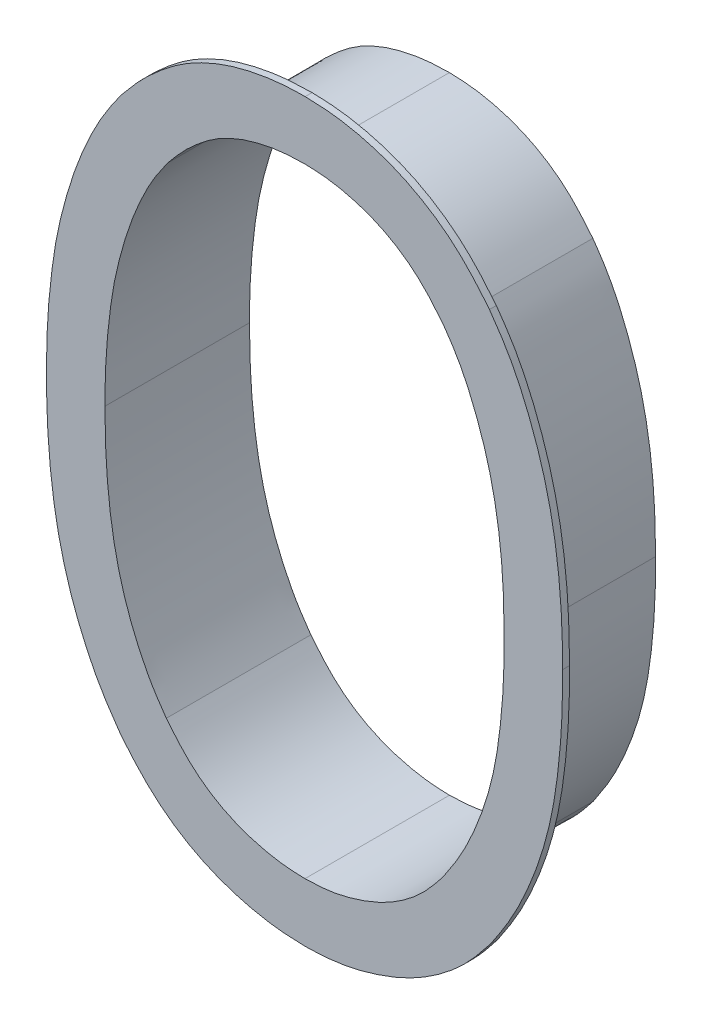
SolidWorks part; units mm, degrees
ref_plane "Front Plane" through (0, 0, 0) normal (0, 0, 1) x (1, 0, 0)
ref_plane "Top Plane" through (0, 0, 0) normal (0, 1, 0) x (1, 0, 0)
ref_plane "Right Plane" through (0, 0, 0) normal (1, 0, 0) x (0, 0, -1)
sketch "Sketch1" plane through (0, 0, 0) normal (0, 0, 1) x (1, 0, 0)
  spline S44 degree 3 poles (5623.5923, 1361.6442) (2863.8993, -1686.6739) (2899.6289, -1569.0458) (2864.1682, -1530.1087) (2863.2577, -1529.2047) (2861.3204, -1527.5284) (2860.2917, -1526.7583) (2858.6691, -1525.6932) (2858.1155, -1525.3526) (2856.9825, -1524.7006) (2856.4033, -1524.39) (2853.4876, -1522.9419) (2851.0525, -1522.1041) (2847.9067, -1521.3759) (2847.2726, -1521.2455) (2845.9931, -1521.0204) (2845.3463, -1520.9257) (2844.0448, -1520.7799) (2843.3925, -1520.731) (2799.3471, -1518.3703) (2752.0518, -1577.1712) (2967.2806, 2475.6155) knots -4.859202 -4.859202 -4.859202 -4.859202 0.125 0.125 0.25 0.25 0.375 0.375 0.4375 0.4375 0.5 0.5 0.75 0.75 0.8125 0.8125 0.875 0.875 0.9375 0.9375 5.089551 5.089551 5.089551 5.089551 only from (2867.551, -1534.0183) to (2840.7781, -1520.6183)
  spline S45 degree 3 poles (2247.577, 2433.1947) (2952.4557, -1632.7722) (2883.5094, -1516.3995) (2835.6295, -1520.9169) (2834.3662, -1521.1201) (2831.8611, -1521.6433) (2830.6199, -1521.9667) (2828.1701, -1522.7885) (2826.9533, -1523.2872) (2824.6238, -1524.4171) (2823.5067, -1525.0559) (2821.3834, -1526.5056) (2820.373, -1527.3102) (2818.8979, -1528.5798) (2818.4133, -1529.0159) (2817.4725, -1529.9117) (2817.0159, -1530.3724) (2783.0829, -1566.7568) (2832.1655, -1679.1716) (-214.1206, 1076.2786) knots -4.430772 -4.430772 -4.430772 -4.430772 0.125 0.125 0.25 0.25 0.375 0.375 0.5 0.5 0.625 0.625 0.75 0.75 0.8125 0.8125 0.875 0.875 5.60901 5.60901 5.60901 5.60901 only from (2840.7781, -1520.6183) to (2814.035, -1533.797)
  spline S46 degree 3 poles (-717.5542, 340.1215) (2932.6815, -1487.8387) (2839.4543, -1495.7986) (2812.0173, -1536.7207) (2811.5485, -1537.469) (2810.6725, -1538.9955) (2810.2643, -1539.7732) (2809.4885, -1541.3484) (2809.1198, -1542.1453) (2808.4177, -1543.7564) (2808.0848, -1544.5707) (2807.4575, -1546.2181) (2807.1635, -1547.0514) (2806.6096, -1548.7344) (2806.3492, -1549.5854) (2805.858, -1551.2934) (2805.6265, -1552.1502) (2805.1979, -1553.8711) (2805.0009, -1554.735) (2804.6469, -1556.4711) (2804.4907, -1557.3434) (2804.2115, -1559.0949) (2804.0885, -1559.974) (2803.866, -1561.7371) (2803.7655, -1562.6207) (2803.4981, -1565.2719) (2803.369, -1567.0422) (2800.0394, -1646.5144) (2893.3062, -1729.7043) (-1191.6183, -1575.2053) knots -3.34907 -3.34907 -3.34907 -3.34907 0.0625 0.0625 0.125 0.125 0.1875 0.1875 0.25 0.25 0.3125 0.3125 0.375 0.375 0.4375 0.4375 0.5 0.5 0.5625 0.5625 0.625 0.625 0.6875 0.6875 0.75 0.75 0.875 0.875 6.351779 6.351779 6.351779 6.351779 only from (2814.035, -1533.797) to (2803.1718, -1574.1413)
  spline S47 degree 3 poles (-1190.6479, -1519.1116) (2887.1329, -1411.3146) (2800.1634, -1497.462) (2803.3576, -1581.1698) (2803.4692, -1582.9239) (2803.794, -1586.4274) (2804.003, -1588.1737) (2804.54, -1591.6435) (2804.8713, -1593.3676) (2805.4826, -1595.934) (2805.7053, -1596.7875) (2806.186, -1598.4752) (2806.4442, -1599.3108) (2807.2746, -1601.7917) (2807.9038, -1603.4105) (2808.9555, -1605.7888) (2809.3231, -1606.5736) (2810.0953, -1608.1261) (2810.501, -1608.8933) (2811.3679, -1610.4019) (2811.8304, -1611.1428) (2839.7617, -1653.2512) (2931.4518, -1664.8342) (-749.5731, -3426.131) knots -5.708122 -5.708122 -5.708122 -5.708122 0.125 0.125 0.25 0.25 0.375 0.375 0.5 0.5 0.5625 0.5625 0.625 0.625 0.75 0.75 0.8125 0.8125 0.875 0.875 0.9375 0.9375 4.477312 4.477312 4.477312 4.477312 only from (2803.1718, -1574.1413) to (2813.8078, -1614.047)
  spline S48 degree 3 poles (29.5815, -4482.6192) (2822.6625, -1460.5193) (2782.5191, -1579.7715) (2817.1933, -1617.9946) (2818.1119, -1618.9015) (2820.0579, -1620.5946) (2821.0854, -1621.3806) (2822.714, -1622.4629) (2823.2715, -1622.8074) (2824.4164, -1623.4634) (2824.9978, -1623.7715) (2827.9332, -1625.2119) (2830.3847, -1626.0579) (2833.5582, -1626.7919) (2834.1982, -1626.9227) (2835.4907, -1627.1478) (2836.1444, -1627.2421) (2883.2083, -1632.4329) (2938.7329, -1513.2193) (2684.2688, -5622.4333) knots -4.727596 -4.727596 -4.727596 -4.727596 0.125 0.125 0.25 0.25 0.375 0.375 0.4375 0.4375 0.5 0.5 0.75 0.75 0.8125 0.8125 0.875 0.875 5.309747 5.309747 5.309747 5.309747 only from (2813.8078, -1614.047) to (2840.7375, -1627.5482)
  spline S49 degree 3 poles (3450.4306, -5578.8149) (2728.9569, -1514.3675) (2798.4471, -1632.3654) (2845.9653, -1627.1771) (2847.2467, -1626.9495) (2849.7793, -1626.334) (2851.0306, -1625.9471) (2852.8911, -1625.2792) (2853.5091, -1625.0402) (2854.7211, -1624.5285) (2855.3168, -1624.2552) (2857.0699, -1623.3772) (2858.1949, -1622.7176) (2859.8236, -1621.628) (2860.3565, -1621.2477) (2861.4006, -1620.4504) (2861.9135, -1620.032) (2863.405, -1618.729) (2864.3347, -1617.8006) (2898.0596, -1579.9006) (2847.2007, -1465.7236) (5901.4164, -4217.2551) knots -4.32716 -4.32716 -4.32716 -4.32716 0.125 0.125 0.25 0.25 0.375 0.375 0.4375 0.4375 0.5 0.5 0.625 0.625 0.6875 0.6875 0.75 0.75 0.875 0.875 5.579937 5.579937 5.579937 5.579937 only from (2840.7375, -1627.5482) to (2867.7085, -1613.7687)
  spline S50 degree 3 poles (6410.7456, -3464.8007) (2752.8813, -1673.5541) (2840.2273, -1656.4052) (2869.6305, -1610.8521) (2870.0866, -1610.1113) (2871.3803, -1607.8538) (2872.151, -1606.3053) (2873.5516, -1603.1417) (2874.1815, -1601.5265) (2875.02, -1599.0533) (2875.2815, -1598.2204) (2875.7661, -1596.5364) (2875.9885, -1595.6886) (2876.594, -1593.137) (2876.9133, -1591.4206) (2877.297, -1588.8288) (2877.4093, -1587.962) (2877.6122, -1586.2245) (2877.7035, -1585.3535) (2877.9422, -1582.7399) (2878.0517, -1580.9952) (2880.8027, -1499.4274) (2790.3135, -1415.3217) (6872.3495, -1523.0841) knots -3.760505 -3.760505 -3.760505 -3.760505 0.0625 0.0625 0.125 0.125 0.25 0.25 0.375 0.375 0.4375 0.4375 0.5 0.5 0.625 0.625 0.6875 0.6875 0.75 0.75 0.875 0.875 6.586269 6.586269 6.586269 6.586269 only from (2867.7085, -1613.7687) to (2878.1982, -1574.0031)
  spline S51 degree 3 poles (6872.2063, -1616.6851) (2793.1681, -1735.7776) (2881.3055, -1650.0072) (2878.0038, -1566.9717) (2877.8888, -1565.2172) (2877.5502, -1561.7134) (2877.3294, -1559.9672) (2876.7655, -1556.5002) (2876.4225, -1554.7778) (2875.8011, -1552.2135) (2875.5756, -1551.3605) (2875.0889, -1549.6722) (2874.8279, -1548.8362) (2873.9969, -1546.3501) (2873.3834, -1544.7202) (2872.3627, -1542.3215) (2872.0054, -1541.5298) (2871.2487, -1539.9657) (2870.8489, -1539.1936) (2869.9897, -1537.6767) (2869.5292, -1536.9325) (2842.2715, -1495.6479) (2749.9543, -1485.2621) (6437.7085, 264.8424) knots -5.658153 -5.658153 -5.658153 -5.658153 0.125 0.125 0.25 0.25 0.375 0.375 0.5 0.5 0.5625 0.5625 0.625 0.625 0.75 0.75 0.8125 0.8125 0.875 0.875 0.9375 0.9375 4.393613 4.393613 4.393613 4.393613 only from (2878.1982, -1574.0031) to (2867.551, -1534.0183)
  spline S52 degree 3 poles (2867.551, -1534.0183) (2866.7267, -1533.0167) (2865.9033, -1532.014) (2864.1682, -1530.1087) (2863.2577, -1529.2047) (2861.3204, -1527.5284) (2860.2917, -1526.7583) (2858.6691, -1525.6932) (2858.1155, -1525.3526) (2856.9825, -1524.7006) (2856.4033, -1524.39) (2853.4876, -1522.9419) (2851.0525, -1522.1041) (2847.9067, -1521.3759) (2847.2726, -1521.2455) (2845.9931, -1521.0204) (2845.3463, -1520.9257) (2844.0448, -1520.7799) (2843.3925, -1520.731) (2842.0862, -1520.661) (2841.4321, -1520.6398) (2840.7781, -1520.6183) knots 0 0 0 0 0.125 0.125 0.25 0.25 0.375 0.375 0.4375 0.4375 0.5 0.5 0.75 0.75 0.8125 0.8125 0.875 0.875 0.9375 0.9375 1 1 1 1
  spline S53 degree 3 poles (2840.7781, -1520.6183) (2839.4823, -1520.646) (2838.1868, -1520.6757) (2835.6295, -1520.9169) (2834.3662, -1521.1201) (2831.8611, -1521.6433) (2830.6199, -1521.9667) (2828.1701, -1522.7885) (2826.9533, -1523.2872) (2824.6238, -1524.4171) (2823.5067, -1525.0559) (2821.3834, -1526.5056) (2820.373, -1527.3102) (2818.8979, -1528.5798) (2818.4133, -1529.0159) (2817.4725, -1529.9117) (2817.0159, -1530.3724) (2815.6894, -1531.7947) (2814.8627, -1532.7963) (2814.035, -1533.797) knots 0 0 0 0 0.125 0.125 0.25 0.25 0.375 0.375 0.5 0.5 0.625 0.625 0.75 0.75 0.8125 0.8125 0.875 0.875 1 1 1 1
  spline S54 degree 3 poles (2814.035, -1533.797) (2813.5203, -1534.5229) (2813.0045, -1535.2483) (2812.0173, -1536.7207) (2811.5485, -1537.469) (2810.6725, -1538.9955) (2810.2643, -1539.7732) (2809.4885, -1541.3484) (2809.1198, -1542.1453) (2808.4177, -1543.7564) (2808.0848, -1544.5707) (2807.4575, -1546.2181) (2807.1635, -1547.0514) (2806.6096, -1548.7344) (2806.3492, -1549.5854) (2805.858, -1551.2934) (2805.6265, -1552.1502) (2805.1979, -1553.8711) (2805.0009, -1554.735) (2804.6469, -1556.4711) (2804.4907, -1557.3434) (2804.2115, -1559.0949) (2804.0885, -1559.974) (2803.866, -1561.7371) (2803.7655, -1562.6207) (2803.4981, -1565.2719) (2803.369, -1567.0422) (2803.2204, -1570.5889) (2803.1964, -1572.3651) (2803.1718, -1574.1413) knots 0 0 0 0 0.0625 0.0625 0.125 0.125 0.1875 0.1875 0.25 0.25 0.3125 0.3125 0.375 0.375 0.4375 0.4375 0.5 0.5 0.5625 0.5625 0.625 0.625 0.6875 0.6875 0.75 0.75 0.875 0.875 1 1 1 1
  spline S55 degree 3 poles (2803.1718, -1574.1413) (2803.1979, -1575.8994) (2803.2236, -1577.6575) (2803.3576, -1581.1698) (2803.4692, -1582.9239) (2803.794, -1586.4274) (2804.003, -1588.1737) (2804.54, -1591.6435) (2804.8713, -1593.3676) (2805.4826, -1595.934) (2805.7053, -1596.7875) (2806.186, -1598.4752) (2806.4442, -1599.3108) (2807.2746, -1601.7917) (2807.9038, -1603.4105) (2808.9555, -1605.7888) (2809.3231, -1606.5736) (2810.0953, -1608.1261) (2810.501, -1608.8933) (2811.3679, -1610.4019) (2811.8304, -1611.1428) (2812.7996, -1612.6039) (2813.3043, -1613.3252) (2813.8078, -1614.047) knots 0 0 0 0 0.125 0.125 0.25 0.25 0.375 0.375 0.5 0.5 0.5625 0.5625 0.625 0.625 0.75 0.75 0.8125 0.8125 0.875 0.875 0.9375 0.9375 1 1 1 1
  spline S56 degree 3 poles (2813.8078, -1614.047) (2814.6301, -1615.0606) (2815.4518, -1616.0749) (2817.1933, -1617.9946) (2818.1119, -1618.9015) (2820.0579, -1620.5946) (2821.0854, -1621.3806) (2822.714, -1622.4629) (2823.2715, -1622.8074) (2824.4164, -1623.4634) (2824.9978, -1623.7715) (2827.9332, -1625.2119) (2830.3847, -1626.0579) (2833.5582, -1626.7919) (2834.1982, -1626.9227) (2835.4907, -1627.1478) (2836.1444, -1627.2421) (2838.1066, -1627.4585) (2839.422, -1627.504) (2840.7375, -1627.5482) knots 0 0 0 0 0.125 0.125 0.25 0.25 0.375 0.375 0.4375 0.4375 0.5 0.5 0.75 0.75 0.8125 0.8125 0.875 0.875 1 1 1 1
  spline S57 degree 3 poles (2840.7375, -1627.5482) (2842.0538, -1627.5052) (2843.3699, -1627.4605) (2845.9653, -1627.1771) (2847.2467, -1626.9495) (2849.7793, -1626.334) (2851.0306, -1625.9471) (2852.8911, -1625.2792) (2853.5091, -1625.0402) (2854.7211, -1624.5285) (2855.3168, -1624.2552) (2857.0699, -1623.3772) (2858.1949, -1622.7176) (2859.8236, -1621.628) (2860.3565, -1621.2477) (2861.4006, -1620.4504) (2861.9135, -1620.032) (2863.405, -1618.729) (2864.3347, -1617.8006) (2866.0803, -1615.8389) (2866.894, -1614.8035) (2867.7085, -1613.7687) knots 0 0 0 0 0.125 0.125 0.25 0.25 0.375 0.375 0.4375 0.4375 0.5 0.5 0.625 0.625 0.6875 0.6875 0.75 0.75 0.875 0.875 1 1 1 1
  spline S58 degree 3 poles (2867.7085, -1613.7687) (2868.196, -1613.0429) (2868.6846, -1612.3176) (2869.6305, -1610.8521) (2870.0866, -1610.1113) (2871.3803, -1607.8538) (2872.151, -1606.3053) (2873.5516, -1603.1417) (2874.1815, -1601.5265) (2875.02, -1599.0533) (2875.2815, -1598.2204) (2875.7661, -1596.5364) (2875.9885, -1595.6886) (2876.594, -1593.137) (2876.9133, -1591.4206) (2877.297, -1588.8288) (2877.4093, -1587.962) (2877.6122, -1586.2245) (2877.7035, -1585.3535) (2877.9422, -1582.7399) (2878.0517, -1580.9952) (2878.1695, -1577.5012) (2878.1838, -1575.7522) (2878.1982, -1574.0031) knots 0 0 0 0 0.0625 0.0625 0.125 0.125 0.25 0.25 0.375 0.375 0.4375 0.4375 0.5 0.5 0.625 0.625 0.6875 0.6875 0.75 0.75 0.875 0.875 1 1 1 1
  spline S59 degree 3 poles (2878.1982, -1574.0031) (2878.1707, -1572.2442) (2878.1435, -1570.4853) (2878.0038, -1566.9717) (2877.8888, -1565.2172) (2877.5502, -1561.7134) (2877.3294, -1559.9672) (2876.7655, -1556.5002) (2876.4225, -1554.7778) (2875.8011, -1552.2135) (2875.5756, -1551.3605) (2875.0889, -1549.6722) (2874.8279, -1548.8362) (2873.9969, -1546.3501) (2873.3834, -1544.7202) (2872.3627, -1542.3215) (2872.0054, -1541.5298) (2871.2487, -1539.9657) (2870.8489, -1539.1936) (2869.9897, -1537.6767) (2869.5292, -1536.9325) (2868.5609, -1535.4658) (2868.0553, -1534.7423) (2867.551, -1534.0183) knots 0 0 0 0 0.125 0.125 0.25 0.25 0.375 0.375 0.5 0.5 0.5625 0.5625 0.625 0.625 0.75 0.75 0.8125 0.8125 0.875 0.875 0.9375 0.9375 1 1 1 1
  spline S60 degree 3 poles (5660.2756, 1313.3797) (2856.4156, -1670.0709) (2887.4383, -1571.0474) (2857.1997, -1537.2991) (2856.5657, -1536.6519) (2855.2096, -1535.4534) (2854.483, -1534.907) (2853.333, -1534.1526) (2852.9388, -1533.9105) (2852.1386, -1533.4513) (2851.7339, -1533.2351) (2849.6859, -1532.2244) (2847.967, -1531.6483) (2845.7445, -1531.1415) (2845.2965, -1531.0503) (2844.3916, -1530.8934) (2843.9341, -1530.8276) (2807.0392, -1526.9137) (2762.8326, -1629.8973) (3023.7967, 2463.9175) knots -5.981424 -5.981424 -5.981424 -5.981424 0.125 0.125 0.25 0.25 0.375 0.375 0.4375 0.4375 0.5 0.5 0.75 0.75 0.8125 0.8125 0.875 0.875 5.850323 5.850323 5.850323 5.850323 only from (2859.5746, -1540.0629) to (2840.7203, -1530.6218)
  spline S61 degree 3 poles (2190.3612, 2414.788) (2932.4724, -1625.4573) (2875.4674, -1527.5067) (2837.1026, -1530.8157) (2836.2158, -1530.9557) (2834.4571, -1531.3119) (2833.5851, -1531.5283) (2832.2956, -1531.9489) (2831.8689, -1532.105) (2831.0212, -1532.4472) (2830.599, -1532.6341) (2829.7754, -1533.0317) (2829.3725, -1533.2435) (2828.5898, -1533.7002) (2828.2106, -1533.9462) (2827.4736, -1534.469) (2827.115, -1534.7447) (2826.4092, -1535.3125) (2826.0618, -1535.6045) (2825.3772, -1536.2028) (2825.0398, -1536.5106) (2824.3831, -1537.1453) (2824.0649, -1537.4718) (2795.8206, -1568.2501) (2838.5799, -1662.5578) (-224.8764, 1049.2327) knots -5.08552 -5.08552 -5.08552 -5.08552 0.125 0.125 0.25 0.25 0.375 0.375 0.4375 0.4375 0.5 0.5 0.5625 0.5625 0.625 0.625 0.6875 0.6875 0.75 0.75 0.8125 0.8125 0.875 0.875 6.543198 6.543198 6.543198 6.543198 only from (2840.7203, -1530.6218) to (2821.9777, -1539.8839)
  spline S62 degree 3 poles (-727.4015, 300.4209) (2936.1542, -1504.8438) (2843.8573, -1506.6945) (2820.2791, -1542.3654) (2819.8914, -1543.0036) (2819.1758, -1544.3086) (2818.8435, -1544.9733) (2818.209, -1546.3172) (2817.9075, -1546.9967) (2817.3363, -1548.371) (2817.0671, -1549.0661) (2816.5625, -1550.4723) (2816.3264, -1551.1833) (2815.8805, -1552.6177) (2815.6704, -1553.3406) (2815.2741, -1554.789) (2815.0885, -1555.5158) (2814.7486, -1556.9755) (2814.5945, -1557.7086) (2814.3216, -1559.182) (2814.0818, -1560.662) (2813.8902, -1562.1517) (2813.7142, -1563.6447) (2813.6344, -1564.392) (2813.4246, -1566.6349) (2813.326, -1568.1325) (2810.506, -1643.9918) (2893.5388, -1723.0667) (-1182.0259, -1573.5803) knots -3.438098 -3.438098 -3.438098 -3.438098 0.0625 0.0625 0.125 0.125 0.1875 0.1875 0.25 0.25 0.3125 0.3125 0.375 0.375 0.4375 0.4375 0.5 0.5 0.5625 0.5625 0.625 0.6875 0.6875 0.75 0.75 0.875 0.875 7.071853 7.071853 7.071853 7.071853 only from (2821.9777, -1539.8839) to (2813.1728, -1574.1361)
  spline S63 degree 3 poles (-1181.2706, -1546.3912) (2887.675, -1416.5356) (2810.5862, -1499.6135) (2813.318, -1580.0797) (2813.4015, -1581.5631) (2813.6509, -1584.5258) (2813.8134, -1586.0068) (2814.2282, -1588.9495) (2814.4829, -1590.412) (2814.9602, -1592.588) (2815.135, -1593.3104) (2815.5169, -1594.7491) (2815.7241, -1595.4649) (2816.3921, -1597.5859) (2816.9027, -1598.9692) (2817.7651, -1600.9987) (2818.0681, -1601.6679) (2818.7041, -1602.9921) (2819.0369, -1603.6473) (2819.7507, -1604.9348) (2820.1357, -1605.5654) (2844.5896, -1642.8286) (2934.6392, -1648.3837) (-738.7814, -3426.5624) knots -6.522514 -6.522514 -6.522514 -6.522514 0.125 0.125 0.25 0.25 0.375 0.375 0.5 0.5 0.5625 0.5625 0.625 0.625 0.75 0.75 0.8125 0.8125 0.875 0.875 0.9375 0.9375 4.630211 4.630211 4.630211 4.630211 only from (2813.1728, -1574.1361) to (2821.8019, -1608.0282)
  spline S64 degree 3 poles (59.4659, -4498.658) (2828.2394, -1477.1161) (2794.9991, -1578.0624) (2824.1716, -1610.8143) (2824.8097, -1611.4599) (2826.1645, -1612.6635) (2826.8816, -1613.2211) (2828.0219, -1613.9855) (2828.4129, -1614.2281) (2829.217, -1614.6888) (2829.63, -1614.9068) (2831.7079, -1615.9191) (2833.4418, -1616.5047) (2835.6792, -1617.0174) (2836.1301, -1617.1091) (2837.0403, -1617.2667) (2837.5008, -1617.3326) (2874.8062, -1621.3093) (2918.7941, -1517.9055) (2683.3129, -5613.0295) knots -5.762777 -5.762777 -5.762777 -5.762777 0.125 0.125 0.25 0.25 0.375 0.375 0.4375 0.4375 0.5 0.5 0.75 0.75 0.8125 0.8125 0.875 0.875 5.861842 5.861842 5.861842 5.861842 only from (2821.8019, -1608.0282) to (2840.7421, -1617.5427)
  spline S65 degree 3 poles (3581.9916, -5546.8161) (2747.4521, -1520.0572) (2806.8426, -1621.216) (2844.4064, -1617.292) (2845.3015, -1617.1326) (2847.0672, -1616.7005) (2847.9381, -1616.4294) (2849.2329, -1615.9689) (2849.6623, -1615.8057) (2850.5154, -1615.4522) (2850.9397, -1615.261) (2852.1792, -1614.6466) (2852.9693, -1614.1827) (2854.4891, -1613.1648) (2855.2177, -1612.6091) (2856.2554, -1611.6929) (2856.5931, -1611.3732) (2857.2446, -1610.7152) (2857.559, -1610.3764) (2885.1835, -1578.8353) (2839.8476, -1484.1867) (5949.7664, -4145.2243) knots -4.915114 -4.915114 -4.915114 -4.915114 0.125 0.125 0.25 0.25 0.375 0.375 0.4375 0.4375 0.5 0.5 0.625 0.625 0.75 0.75 0.8125 0.8125 0.875 0.875 6.483637 6.483637 6.483637 6.483637 only from (2840.7421, -1617.5427) to (2859.6176, -1607.8798)
  spline S66 degree 3 poles (6296.3594, -3650.1271) (2750.3486, -1655.8584) (2834.6811, -1646.8437) (2861.2472, -1605.3955) (2861.6324, -1604.7624) (2862.719, -1602.825) (2863.3633, -1601.4896) (2864.2407, -1599.4379) (2864.5177, -1598.7455) (2865.0366, -1597.356) (2865.2795, -1596.6574) (2865.9568, -1594.5497) (2866.3386, -1593.1284) (2866.9634, -1590.2539) (2867.206, -1588.8005) (2867.5009, -1586.6044) (2867.5885, -1585.8699) (2867.7482, -1584.3973) (2867.8198, -1583.6588) (2867.9434, -1582.1818) (2867.9957, -1581.4428) (2868.0781, -1579.9641) (2868.108, -1579.2242) (2870.3618, -1502.3714) (2790.1224, -1422.7773) (6862.7887, -1518.4977) knots -4.020864 -4.020864 -4.020864 -4.020864 0.0625 0.0625 0.125 0.125 0.25 0.25 0.3125 0.3125 0.375 0.375 0.5 0.5 0.625 0.625 0.6875 0.6875 0.75 0.75 0.8125 0.8125 0.875 0.875 7.301658 7.301658 7.301658 7.301658 only from (2859.6176, -1607.8798) to (2868.1976, -1574.0402)
  spline S67 degree 3 poles (6862.87, -1587.6778) (2793.0545, -1730.2157) (2870.8559, -1647.7121) (2868.0461, -1568.0938) (2867.9601, -1566.6098) (2867.7007, -1563.6466) (2867.5297, -1562.1653) (2867.0912, -1559.2241) (2866.8232, -1557.7631) (2866.3344, -1555.5888) (2866.157, -1554.8669) (2865.7702, -1553.4293) (2865.5601, -1552.7133) (2864.8877, -1550.589) (2864.3858, -1549.1977) (2863.5542, -1547.1474) (2863.263, -1546.4705) (2862.6467, -1545.1325) (2862.322, -1544.4712) (2861.6208, -1543.1727) (2861.2399, -1542.5376) (2837.7601, -1506.4357) (2745.8952, -1502.9761) (6430.4921, 258.2368) knots -6.448256 -6.448256 -6.448256 -6.448256 0.125 0.125 0.25 0.25 0.375 0.375 0.5 0.5 0.5625 0.5625 0.625 0.625 0.75 0.75 0.8125 0.8125 0.875 0.875 0.9375 0.9375 4.493008 4.493008 4.493008 4.493008 only from (2868.1976, -1574.0402) to (2859.5746, -1540.0629)
  spline S68 degree 3 poles (2859.5746, -1540.0629) (2858.994, -1539.3577) (2858.4128, -1538.6531) (2857.1997, -1537.2991) (2856.5657, -1536.6519) (2855.2096, -1535.4534) (2854.483, -1534.907) (2853.333, -1534.1526) (2852.9388, -1533.9105) (2852.1386, -1533.4513) (2851.7339, -1533.2351) (2849.6859, -1532.2244) (2847.967, -1531.6483) (2845.7445, -1531.1415) (2845.2965, -1531.0503) (2844.3916, -1530.8934) (2843.9341, -1530.8276) (2842.5609, -1530.6819) (2841.6405, -1530.6523) (2840.7203, -1530.6218) knots 0 0 0 0 0.125 0.125 0.25 0.25 0.375 0.375 0.4375 0.4375 0.5 0.5 0.75 0.75 0.8125 0.8125 0.875 0.875 1 1 1 1
  spline S69 degree 3 poles (2840.7203, -1530.6218) (2839.8103, -1530.6414) (2838.9002, -1530.6607) (2837.1026, -1530.8157) (2836.2158, -1530.9557) (2834.4571, -1531.3119) (2833.5851, -1531.5283) (2832.2956, -1531.9489) (2831.8689, -1532.105) (2831.0212, -1532.4472) (2830.599, -1532.6341) (2829.7754, -1533.0317) (2829.3725, -1533.2435) (2828.5898, -1533.7002) (2828.2106, -1533.9462) (2827.4736, -1534.469) (2827.115, -1534.7447) (2826.4092, -1535.3125) (2826.0618, -1535.6045) (2825.3772, -1536.2028) (2825.0398, -1536.5106) (2824.3831, -1537.1453) (2824.0649, -1537.4718) (2823.1408, -1538.4788) (2822.5591, -1539.1812) (2821.9777, -1539.8839) knots 0 0 0 0 0.125 0.125 0.25 0.25 0.375 0.375 0.4375 0.4375 0.5 0.5 0.5625 0.5625 0.625 0.625 0.6875 0.6875 0.75 0.75 0.8125 0.8125 0.875 0.875 1 1 1 1
  spline S70 degree 3 poles (2821.9777, -1539.8839) (2821.5418, -1540.4989) (2821.1062, -1541.114) (2820.2791, -1542.3654) (2819.8914, -1543.0036) (2819.1758, -1544.3086) (2818.8435, -1544.9733) (2818.209, -1546.3172) (2817.9075, -1546.9967) (2817.3363, -1548.371) (2817.0671, -1549.0661) (2816.5625, -1550.4723) (2816.3264, -1551.1833) (2815.8805, -1552.6177) (2815.6704, -1553.3406) (2815.2741, -1554.789) (2815.0885, -1555.5158) (2814.7486, -1556.9755) (2814.5945, -1557.7086) (2814.3216, -1559.182) (2814.0818, -1560.662) (2813.8902, -1562.1517) (2813.7142, -1563.6447) (2813.6344, -1564.392) (2813.4246, -1566.6349) (2813.326, -1568.1325) (2813.2144, -1571.1324) (2813.1936, -1572.6343) (2813.1728, -1574.1361) knots 0 0 0 0 0.0625 0.0625 0.125 0.125 0.1875 0.1875 0.25 0.25 0.3125 0.3125 0.375 0.375 0.4375 0.4375 0.5 0.5 0.5625 0.5625 0.625 0.6875 0.6875 0.75 0.75 0.875 0.875 1 1 1 1
  spline S71 degree 3 poles (2813.1728, -1574.1361) (2813.1949, -1575.6228) (2813.2171, -1577.1094) (2813.318, -1580.0797) (2813.4015, -1581.5631) (2813.6509, -1584.5258) (2813.8134, -1586.0068) (2814.2282, -1588.9495) (2814.4829, -1590.412) (2814.9602, -1592.588) (2815.135, -1593.3104) (2815.5169, -1594.7491) (2815.7241, -1595.4649) (2816.3921, -1597.5859) (2816.9027, -1598.9692) (2817.7651, -1600.9987) (2818.0681, -1601.6679) (2818.7041, -1602.9921) (2819.0369, -1603.6473) (2819.7507, -1604.9348) (2820.1357, -1605.5654) (2820.9497, -1606.8058) (2821.3756, -1607.417) (2821.8019, -1608.0282) knots 0 0 0 0 0.125 0.125 0.25 0.25 0.375 0.375 0.5 0.5 0.5625 0.5625 0.625 0.625 0.75 0.75 0.8125 0.8125 0.875 0.875 0.9375 0.9375 1 1 1 1
  spline S72 degree 3 poles (2821.8019, -1608.0282) (2822.38, -1608.7406) (2822.9586, -1609.4525) (2824.1716, -1610.8143) (2824.8097, -1611.4599) (2826.1645, -1612.6635) (2826.8816, -1613.2211) (2828.0219, -1613.9855) (2828.4129, -1614.2281) (2829.217, -1614.6888) (2829.63, -1614.9068) (2831.7079, -1615.9191) (2833.4418, -1616.5047) (2835.6792, -1617.0174) (2836.1301, -1617.1091) (2837.0403, -1617.2667) (2837.5008, -1617.3326) (2838.8861, -1617.4803) (2839.8141, -1617.5113) (2840.7421, -1617.5427) knots 0 0 0 0 0.125 0.125 0.25 0.25 0.375 0.375 0.4375 0.4375 0.5 0.5 0.75 0.75 0.8125 0.8125 0.875 0.875 1 1 1 1
  spline S73 degree 3 poles (2840.7421, -1617.5427) (2841.6652, -1617.5123) (2842.5882, -1617.4819) (2844.4064, -1617.292) (2845.3015, -1617.1326) (2847.0672, -1616.7005) (2847.9381, -1616.4294) (2849.2329, -1615.9689) (2849.6623, -1615.8057) (2850.5154, -1615.4522) (2850.9397, -1615.261) (2852.1792, -1614.6466) (2852.9693, -1614.1827) (2854.4891, -1613.1648) (2855.2177, -1612.6091) (2856.2554, -1611.6929) (2856.5931, -1611.3732) (2857.2446, -1610.7152) (2857.559, -1610.3764) (2858.4724, -1609.3336) (2859.0452, -1608.6068) (2859.6176, -1607.8798) knots 0 0 0 0 0.125 0.125 0.25 0.25 0.375 0.375 0.4375 0.4375 0.5 0.5 0.625 0.625 0.75 0.75 0.8125 0.8125 0.875 0.875 1 1 1 1
  spline S74 degree 3 poles (2859.6176, -1607.8798) (2860.0321, -1607.2626) (2860.4462, -1606.6452) (2861.2472, -1605.3955) (2861.6324, -1604.7624) (2862.719, -1602.825) (2863.3633, -1601.4896) (2864.2407, -1599.4379) (2864.5177, -1598.7455) (2865.0366, -1597.356) (2865.2795, -1596.6574) (2865.9568, -1594.5497) (2866.3386, -1593.1284) (2866.9634, -1590.2539) (2867.206, -1588.8005) (2867.5009, -1586.6044) (2867.5885, -1585.8699) (2867.7482, -1584.3973) (2867.8198, -1583.6588) (2867.9434, -1582.1818) (2867.9957, -1581.4428) (2868.0781, -1579.9641) (2868.108, -1579.2242) (2868.1732, -1577.0036) (2868.1854, -1575.5219) (2868.1976, -1574.0402) knots 0 0 0 0 0.0625 0.0625 0.125 0.125 0.25 0.25 0.3125 0.3125 0.375 0.375 0.5 0.5 0.625 0.625 0.6875 0.6875 0.75 0.75 0.8125 0.8125 0.875 0.875 1 1 1 1
  spline S75 degree 3 poles (2868.1976, -1574.0402) (2868.1743, -1572.5528) (2868.151, -1571.0654) (2868.0461, -1568.0938) (2867.9601, -1566.6098) (2867.7007, -1563.6466) (2867.5297, -1562.1653) (2867.0912, -1559.2241) (2866.8232, -1557.7631) (2866.3344, -1555.5888) (2866.157, -1554.8669) (2865.7702, -1553.4293) (2865.5601, -1552.7133) (2864.8877, -1550.589) (2864.3858, -1549.1977) (2863.5542, -1547.1474) (2863.263, -1546.4705) (2862.6467, -1545.1325) (2862.322, -1544.4712) (2861.6208, -1543.1727) (2861.2399, -1542.5376) (2860.4286, -1541.2903) (2860.0018, -1540.6765) (2859.5746, -1540.0629) knots 0 0 0 0 0.125 0.125 0.25 0.25 0.375 0.375 0.5 0.5 0.5625 0.5625 0.625 0.625 0.75 0.75 0.8125 0.8125 0.875 0.875 0.9375 0.9375 1 1 1 1
  dimension "D1" = 5
  dimension "D2" = 5
extrude "Boss-Extrude1" add sketch "Sketch1" along normal blind 1 and the other way blind 20
sketch3d "3DSketch1"
  spline S0 degree 5 poles (2777.4956, -3616.8164, 1) (2771.5169, -2410.8399, 1) (2779.4982, -1811.9825, 1) (2796.9834, -1616.2173, 1) (2819.4505, -1619.8557, 1) (2841.8118, -1619.0055, 1) (2842.0923, -1618.9932, 1) (2842.7784, -1618.9571, 1) (2843.4636, -1618.9006, 1) (2843.8681, -1618.8589, 1) (2844.7178, -1618.7516, 1) (2845.5605, -1618.5981, 1) (2846.001, -1618.5057, 1) (2846.948, -1618.2826, 1) (2847.8826, -1618.0137, 1) (2848.3813, -1617.8572, 1) (2849.4328, -1617.5018, 1) (2850.4692, -1617.1028, 1) (2851.0114, -1616.8773, 1) (2852.0701, -1616.3978, 1) (2853.0924, -1615.844, 1) (2853.5893, -1615.553, 1) (2854.5058, -1614.977, 1) (2855.3887, -1614.3511, 1) (2855.7938, -1614.047, 1) (2856.5402, -1613.4525, 1) (2857.2519, -1612.8171, 1) (2857.5781, -1612.5103, 1) (2858.1954, -1611.8993, 1) (2858.7821, -1611.2592, 1) (2859.0602, -1610.9434, 1) (2859.5238, -1610.3985, 1) (2859.9747, -1609.8435, 1) (2860.1587, -1609.6136, 1) (2875.759, -1589.9578, 1) (2888.13, -1567.7626, 1) (3057.068, -1669.0583, 1) (3542.583, -2019.2963, 1) (4505.2564, -2743.6565, 1) knots -4.68935 -4.68935 -4.68935 -4.68935 -4.68935 -4.68935 0.021729 0.021729 0.021729 0.081586 0.081586 0.081586 0.168224 0.168224 0.168224 0.264114 0.264114 0.264114 0.375486 0.375486 0.375486 0.500556 0.500556 0.500556 0.623143 0.623143 0.623143 0.731014 0.731014 0.731014 0.826417 0.826417 0.826417 0.91609 0.91609 0.91609 0.978877 0.978877 0.978877 6.266542 6.266542 6.266542 6.266542 6.266542 6.266542 only from (2840.7414, -1619.0435, 1) to (2860.8312, -1608.7631, 1)
  spline S1 degree 5 poles (4397.2962, -2886.5859, 1) (3436.5593, -2157.5568, 1) (2968.1974, -1785.2284, 1) (2826.7415, -1649.5286, 1) (2846.741, -1630.1103, 1) (2861.8868, -1607.1786, 1) (2862.1459, -1606.7792, 1) (2862.7812, -1605.7732, 1) (2863.3742, -1604.7411, 1) (2863.7153, -1604.1135, 1) (2864.3618, -1602.8588, 1) (2864.9561, -1601.5791, 1) (2865.2375, -1600.9415, 1) (2865.783, -1599.6421, 1) (2866.2833, -1598.3247, 1) (2866.5243, -1597.6544, 1) (2866.9814, -1596.3061, 1) (2867.3883, -1594.9416, 1) (2867.5788, -1594.256, 1) (2867.9376, -1592.8622, 1) (2868.2415, -1591.4554, 1) (2868.382, -1590.7413, 1) (2868.6418, -1589.2906, 1) (2868.855, -1587.8327, 1) (2868.9528, -1587.0932, 1) (2869.1331, -1585.5989, 1) (2869.2862, -1584.1016, 1) (2869.3558, -1583.3457, 1) (2869.4795, -1581.8112, 1) (2869.5648, -1580.2739, 1) (2869.5992, -1579.4941, 1) (2869.6433, -1578.189, 1) (2869.6679, -1576.8836, 1) (2869.6754, -1576.3585, 1) (2870.1198, -1537.0073, 1) (2866.1336, -1497.6324, 1) (3060.8935, -1459.8449, 1) (3657.3537, -1424.2043, 1) (4858.0646, -1391.8498, 1) knots -3.675995 -3.675995 -3.675995 -3.675995 -3.675995 -3.675995 0.026102 0.026102 0.026102 0.091367 0.091367 0.091367 0.189244 0.189244 0.189244 0.284775 0.284775 0.284775 0.382411 0.382411 0.382411 0.479937 0.479937 0.479937 0.57969 0.57969 0.57969 0.681959 0.681959 0.681959 0.786036 0.786036 0.786036 0.893054 0.893054 0.893054 0.965071 0.965071 0.965071 6.289432 6.289432 6.289432 6.289432 6.289432 6.289432 only from (2860.8312, -1608.7631, 1) to (2869.6977, -1574.0346, 1)
  spline S2 degree 5 poles (4858.1254, -1755.0559, 1) (3655.9441, -1723.957, 1) (3059.7382, -1688.7669, 1) (2865.8062, -1650.8714, 1) (2870.4516, -1610.9827, 1) (2869.6464, -1571.1306, 1) (2869.6303, -1570.4731, 1) (2869.5796, -1568.8351, 1) (2869.4945, -1567.1982, 1) (2869.4301, -1566.219, 1) (2869.2756, -1564.3013, 1) (2869.0619, -1562.3892, 1) (2868.9423, -1561.4541, 1) (2868.6889, -1559.7051, 1) (2868.3786, -1557.9651, 1) (2868.2206, -1557.1557, 1) (2867.9008, -1555.659, 1) (2867.5288, -1554.1745, 1) (2867.3461, -1553.4926, 1) (2866.9858, -1552.2307, 1) (2866.5871, -1550.9805, 1) (2866.3949, -1550.4053, 1) (2865.9962, -1549.2625, 1) (2865.5683, -1548.1303, 1) (2865.3475, -1547.5682, 1) (2864.9029, -1546.4796, 1) (2864.4297, -1545.4029, 1) (2864.1913, -1544.883, 1) (2863.6903, -1543.8433, 1) (2863.1432, -1542.8265, 1) (2862.8553, -1542.3202, 1) (2862.3577, -1541.4927, 1) (2861.826, -1540.6873, 1) (2861.6112, -1540.3701, 1) (2846.4484, -1518.3361, 1) (2827.3054, -1499.357, 1) (2966.1332, -1359.6153, 1) (3424.2221, -974.8368, 1) (4362.7688, -220.909, 1) knots -5.313434 -5.313434 -5.313434 -5.313434 -5.313434 -5.313434 0.043429 0.043429 0.043429 0.133304 0.133304 0.133304 0.267366 0.267366 0.267366 0.396147 0.396147 0.396147 0.508784 0.508784 0.508784 0.605224 0.605224 0.605224 0.68807 0.68807 0.68807 0.770592 0.770592 0.770592 0.84872 0.84872 0.84872 0.928258 0.928258 0.928258 0.980589 0.980589 0.980589 4.58232 4.58232 4.58232 4.58232 4.58232 4.58232 only from (2869.6977, -1574.0346, 1) to (2860.771, -1539.1562, 1)
  spline S3 degree 5 poles (4483.8943, -373.6882, 1) (3537.3672, -1119.0074, 1) (3058.867, -1478.0491, 1) (2891.1, -1581.7983, 1) (2877.0849, -1558.8399, 1) (2860.0889, -1538.3306, 1) (2859.8978, -1538.1017, 1) (2859.4346, -1537.5532, 1) (2858.9612, -1537.0132, 1) (2858.68, -1536.7014, 1) (2858.094, -1536.0739, 1) (2857.4817, -1535.4716, 1) (2857.1615, -1535.1714, 1) (2856.4622, -1534.5502, 1) (2855.7252, -1533.9737, 1) (2855.3245, -1533.6795, 1) (2854.4547, -1533.0775, 1) (2853.554, -1532.5234, 1) (2853.0682, -1532.2439, 1) (2852.0658, -1531.7065, 1) (2851.0315, -1531.2326, 1) (2850.4994, -1531.0086, 1) (2849.4772, -1530.6149, 1) (2848.4345, -1530.281, 1) (2847.9373, -1530.1355, 1) (2846.9976, -1529.8839, 1) (2846.0488, -1529.6695, 1) (2845.6035, -1529.5786, 1) (2844.7512, -1529.425, 1) (2843.8924, -1529.3131, 1) (2843.4831, -1529.2689, 1) (2842.7963, -1529.2092, 1) (2842.1083, -1529.1724, 1) (2841.831, -1529.1603, 1) (2818.9582, -1528.2961, 1) (2796.0518, -1531.7396, 1) (2774.9738, -1335.8369, 1) (2757.0281, -737.1203, 1) (2744.2626, 467.3929, 1) knots -5.638201 -5.638201 -5.638201 -5.638201 -5.638201 -5.638201 0.020394 0.020394 0.020394 0.084454 0.084454 0.084454 0.174634 0.174634 0.174634 0.268859 0.268859 0.268859 0.375482 0.375482 0.375482 0.495778 0.495778 0.495778 0.619637 0.619637 0.619637 0.730851 0.730851 0.730851 0.828455 0.828455 0.828455 0.916841 0.916841 0.916841 0.97647 0.97647 0.97647 5.833814 5.833814 5.833814 5.833814 5.833814 5.833814 only from (2860.771, -1539.1562, 1) to (2840.729, -1529.1213, 1)
  spline S4 degree 5 poles (2937.7952, 467.2814, 1) (2924.3763, -738.1261, 1) (2906.0109, -1336.7023, 1) (2884.948, -1532.3225, 1) (2862.2723, -1528.5502, 1) (2839.6258, -1529.1476, 1) (2839.3494, -1529.1565, 1) (2838.6635, -1529.1844, 1) (2837.9784, -1529.2326, 1) (2837.57, -1529.2693, 1) (2836.7215, -1529.3637, 1) (2835.8786, -1529.4982, 1) (2835.442, -1529.578, 1) (2834.5064, -1529.7681, 1) (2833.5784, -1529.9934, 1) (2833.0848, -1530.1257, 1) (2832.0668, -1530.4287, 1) (2831.07, -1530.7967, 1) (2830.5589, -1531.0048, 1) (2829.5463, -1531.4563, 1) (2828.5648, -1531.9733, 1) (2828.0815, -1532.2503, 1) (2827.1832, -1532.8123, 1) (2826.3329, -1533.4432, 1) (2825.9379, -1533.7549, 1) (2825.1965, -1534.3667, 1) (2824.4722, -1534.9977, 1) (2824.1325, -1535.3041, 1) (2823.4911, -1535.9077, 1) (2822.8802, -1536.5423, 1) (2822.5926, -1536.8534, 1) (2822.1174, -1537.3855, 1) (2821.6548, -1537.928, 1) (2821.4685, -1538.1496, 1) (2805.2038, -1557.6628, 1) (2791.9959, -1579.7573, 1) (2626.5316, -1472.9026, 1) (2153.2699, -1106.1302, 1) (1215.405, -348.8298, 1) knots -4.811181 -4.811181 -4.811181 -4.811181 -4.811181 -4.811181 0.023777 0.023777 0.023777 0.083545 0.083545 0.083545 0.172095 0.172095 0.172095 0.26794 0.26794 0.26794 0.378236 0.378236 0.378236 0.497314 0.497314 0.497314 0.617444 0.617444 0.617444 0.726031 0.726031 0.726031 0.824839 0.824839 0.824839 0.916329 0.916329 0.916329 0.978889 0.978889 0.978889 6.40556 6.40556 6.40556 6.40556 6.40556 6.40556 only from (2840.729, -1529.1213, 1) to (2820.7864, -1538.9708, 1)
  spline S5 degree 5 poles (1336.661, -200.2848, 1) (2264.0965, -973.0372, 1) (2715.9905, -1365.1543, 1) (2852.5253, -1504.8208, 1) (2833.5171, -1520.5724, 1) (2819.7186, -1540.4944, 1) (2819.4557, -1540.8832, 1) (2818.8128, -1541.8705, 1) (2818.2285, -1542.8937, 1) (2817.895, -1543.52, 1) (2817.2608, -1544.7828, 1) (2816.6738, -1546.0672, 1) (2816.3936, -1546.7117, 1) (2815.8462, -1548.0391, 1) (2815.3516, -1549.3871, 1) (2815.1116, -1550.0801, 1) (2814.6533, -1551.4763, 1) (2814.2356, -1552.8848, 1) (2814.0368, -1553.5933, 1) (2813.6571, -1555.0296, 1) (2813.3221, -1556.4773, 1) (2813.1652, -1557.2106, 1) (2812.8754, -1558.6914, 1) (2812.6409, -1560.1817, 1) (2812.5344, -1560.9332, 1) (2812.3384, -1562.4483, 1) (2812.1689, -1563.9662, 1) (2812.0913, -1564.7307, 1) (2811.9511, -1566.2844, 1) (2811.85, -1567.8413, 1) (2811.808, -1568.632, 1) (2811.7524, -1569.9533, 1) (2811.719, -1571.275, 1) (2811.7082, -1571.8054, 1) (2811.0408, -1611.0448, 1) (2814.8766, -1650.3222, 1) (2620.0219, -1687.3954, 1) (2023.5064, -1721.0848, 1) (822.6941, -1749.9001, 1) knots -3.190055 -3.190055 -3.190055 -3.190055 -3.190055 -3.190055 0.024959 0.024959 0.024959 0.088462 0.088462 0.088462 0.18442 0.18442 0.18442 0.279534 0.279534 0.279534 0.378768 0.378768 0.378768 0.478375 0.478375 0.478375 0.579853 0.579853 0.579853 0.682587 0.682587 0.682587 0.786597 0.786597 0.786597 0.893776 0.893776 0.893776 0.965592 0.965592 0.965592 6.206678 6.206678 6.206678 6.206678 6.206678 6.206678 only from (2820.7864, -1538.9708, 1) to (2811.6727, -1574.1369, 1)
  spline S6 degree 5 poles (824.5918, -1380.4562, 1) (2025.7824, -1417.1234, 1) (2621.5542, -1455.6045, 1) (2815.4649, -1495.2578, 1) (2810.94, -1536.1491, 1) (2811.721, -1577.0249, 1) (2811.7364, -1577.6839, 1) (2811.7848, -1579.3185, 1) (2811.8675, -1580.9518, 1) (2811.9295, -1581.9261, 1) (2812.0773, -1583.8401, 1) (2812.278, -1585.7495, 1) (2812.3906, -1586.6863, 1) (2812.6356, -1588.4772, 1) (2812.9413, -1590.2591, 1) (2813.1024, -1591.1083, 1) (2813.4401, -1592.7197, 1) (2813.8404, -1594.3168, 1) (2814.0451, -1595.0719, 1) (2814.4648, -1596.5079, 1) (2814.9397, -1597.9266, 1) (2815.1787, -1598.5991, 1) (2815.6746, -1599.9159, 1) (2816.2188, -1601.2132, 1) (2816.4985, -1601.8476, 1) (2817.0866, -1603.1183, 1) (2817.7208, -1604.3675, 1) (2818.0552, -1604.9905, 1) (2818.6397, -1606.0113, 1) (2819.2776, -1606.9993, 1) (2819.5385, -1607.3897, 1) (2833.7342, -1628.1691, 1) (2852.9969, -1644.9973, 1) (2715.1447, -1783.7514, 1) (2258.9019, -2170.7908, 1) (1322.6816, -2932.0879, 1) knots -5.461291 -5.461291 -5.461291 -5.461291 -5.461291 -5.461291 0.042971 0.042971 0.042971 0.133176 0.133176 0.133176 0.266741 0.266741 0.266741 0.395827 0.395827 0.395827 0.51404 0.51404 0.51404 0.621055 0.621055 0.621055 0.718685 0.718685 0.718685 0.813533 0.813533 0.813533 0.910209 0.910209 0.910209 0.974441 0.974441 0.974441 4.352101 4.352101 4.352101 4.352101 4.352101 4.352101 only from (2811.6727, -1574.1369, 1) to (2820.6028, -1608.931, 1)
  spline S7 degree 5 poles (1195.9153, -2772.8108, 1) (2143.5952, -2030.6622, 1) (2624.1382, -1671.6356, 1) (2791.9478, -1567.5409, 1) (2805.0649, -1589.9296, 1) (2821.2949, -1609.7806, 1) (2821.4825, -1610.0082, 1) (2821.9411, -1610.5574, 1) (2822.4111, -1611.0973, 1) (2822.6922, -1611.4103, 1) (2823.2812, -1612.0421, 1) (2823.8983, -1612.6469, 1) (2824.2223, -1612.9497, 1) (2824.9269, -1613.5768, 1) (2825.6643, -1614.1657, 1) (2826.064, -1614.4665, 1) (2826.933, -1615.0812, 1) (2827.8397, -1615.6389, 1) (2828.3301, -1615.9188, 1) (2829.3408, -1616.4541, 1) (2830.3824, -1616.9257, 1) (2830.9171, -1617.1484, 1) (2831.9479, -1617.5423, 1) (2832.9985, -1617.8786, 1) (2833.5017, -1618.0261, 1) (2834.4504, -1618.2805, 1) (2835.4085, -1618.4963, 1) (2835.857, -1618.5874, 1) (2836.7167, -1618.741, 1) (2837.5829, -1618.8518, 1) (2837.9965, -1618.8955, 1) (2838.6915, -1618.9547, 1) (2839.3876, -1618.9921, 1) (2839.6689, -1619.0046, 1) (2862.5166, -1619.8871, 1) (2885.4319, -1616.3789, 1) (2904.9941, -1812.2471, 1) (2918.3494, -2411.067, 1) (2921.8985, -3616.1663, 1) knots -5.392037 -5.392037 -5.392037 -5.392037 -5.392037 -5.392037 0.021604 0.021604 0.021604 0.084614 0.084614 0.084614 0.174417 0.174417 0.174417 0.269072 0.269072 0.269072 0.375749 0.375749 0.375749 0.496167 0.496167 0.496167 0.619716 0.619716 0.619716 0.731628 0.731628 0.731628 0.829318 0.829318 0.829318 0.918078 0.918078 0.918078 0.978211 0.978211 0.978211 5.801168 5.801168 5.801168 5.801168 5.801168 5.801168 only from (2820.6028, -1608.931, 1) to (2840.7414, -1619.0435, 1)
  spline S8 degree 5 poles (2840.7414, -1619.0435, 1) (2840.8433, -1619.0401, 1) (2840.9451, -1619.0367, 1) (2841.047, -1619.0333, 1) (2841.4294, -1619.02, 1) (2841.8118, -1619.0055, 1) (2842.0923, -1618.9932, 1) (2842.7784, -1618.9571, 1) (2843.4636, -1618.9006, 1) (2843.8681, -1618.8589, 1) (2844.7178, -1618.7516, 1) (2845.5605, -1618.5981, 1) (2846.001, -1618.5057, 1) (2846.948, -1618.2826, 1) (2847.8826, -1618.0137, 1) (2848.3813, -1617.8572, 1) (2849.4328, -1617.5018, 1) (2850.4692, -1617.1028, 1) (2851.0114, -1616.8773, 1) (2852.0701, -1616.3978, 1) (2853.0924, -1615.844, 1) (2853.5893, -1615.553, 1) (2854.5058, -1614.977, 1) (2855.3887, -1614.3511, 1) (2855.7938, -1614.047, 1) (2856.5402, -1613.4525, 1) (2857.2519, -1612.8171, 1) (2857.5781, -1612.5103, 1) (2858.1954, -1611.8993, 1) (2858.7821, -1611.2592, 1) (2859.0602, -1610.9434, 1) (2859.5238, -1610.3985, 1) (2859.9747, -1609.8435, 1) (2860.1587, -1609.6136, 1) (2860.4034, -1609.3054, 1) (2860.6473, -1608.9965, 1) (2860.7086, -1608.9187, 1) (2860.7699, -1608.8409, 1) (2860.8312, -1608.7631, 1) knots 0 0 0 0 0 0 0.021729 0.021729 0.021729 0.081586 0.081586 0.081586 0.168224 0.168224 0.168224 0.264114 0.264114 0.264114 0.375486 0.375486 0.375486 0.500556 0.500556 0.500556 0.623143 0.623143 0.623143 0.731014 0.731014 0.731014 0.826417 0.826417 0.826417 0.91609 0.91609 0.91609 0.978877 0.978877 0.978877 1 1 1 1 1 1
  spline S9 degree 5 poles (2860.8312, -1608.7631, 1) (2860.9373, -1608.6051, 1) (2861.0434, -1608.447, 1) (2861.1493, -1608.2888, 1) (2861.5195, -1607.7347, 1) (2861.8868, -1607.1786, 1) (2862.1459, -1606.7792, 1) (2862.7812, -1605.7732, 1) (2863.3742, -1604.7411, 1) (2863.7153, -1604.1135, 1) (2864.3618, -1602.8588, 1) (2864.9561, -1601.5791, 1) (2865.2375, -1600.9415, 1) (2865.783, -1599.6421, 1) (2866.2833, -1598.3247, 1) (2866.5243, -1597.6544, 1) (2866.9814, -1596.3061, 1) (2867.3883, -1594.9416, 1) (2867.5788, -1594.256, 1) (2867.9376, -1592.8622, 1) (2868.2415, -1591.4554, 1) (2868.382, -1590.7413, 1) (2868.6418, -1589.2906, 1) (2868.855, -1587.8327, 1) (2868.9528, -1587.0932, 1) (2869.1331, -1585.5989, 1) (2869.2862, -1584.1016, 1) (2869.3558, -1583.3457, 1) (2869.4795, -1581.8112, 1) (2869.5648, -1580.2739, 1) (2869.5992, -1579.4941, 1) (2869.6433, -1578.189, 1) (2869.6679, -1576.8836, 1) (2869.6754, -1576.3585, 1) (2869.6842, -1575.5786, 1) (2869.6913, -1574.7987, 1) (2869.6935, -1574.544, 1) (2869.6956, -1574.2893, 1) (2869.6977, -1574.0346, 1) knots 0 0 0 0 0 0 0.026102 0.026102 0.026102 0.091367 0.091367 0.091367 0.189244 0.189244 0.189244 0.284775 0.284775 0.284775 0.382411 0.382411 0.382411 0.479937 0.479937 0.479937 0.57969 0.57969 0.57969 0.681959 0.681959 0.681959 0.786036 0.786036 0.786036 0.893054 0.893054 0.893054 0.965071 0.965071 0.965071 1 1 1 1 1 1
  spline S10 degree 5 poles (2869.6977, -1574.0346, 1) (2869.6927, -1573.7168, 1) (2869.6877, -1573.3991, 1) (2869.6826, -1573.0813, 1) (2869.6661, -1572.1059, 1) (2869.6464, -1571.1306, 1) (2869.6303, -1570.4731, 1) (2869.5796, -1568.8351, 1) (2869.4945, -1567.1982, 1) (2869.4301, -1566.219, 1) (2869.2756, -1564.3013, 1) (2869.0619, -1562.3892, 1) (2868.9423, -1561.4541, 1) (2868.6889, -1559.7051, 1) (2868.3786, -1557.9651, 1) (2868.2206, -1557.1557, 1) (2867.9008, -1555.659, 1) (2867.5288, -1554.1745, 1) (2867.3461, -1553.4926, 1) (2866.9858, -1552.2307, 1) (2866.5871, -1550.9805, 1) (2866.3949, -1550.4053, 1) (2865.9962, -1549.2625, 1) (2865.5683, -1548.1303, 1) (2865.3475, -1547.5682, 1) (2864.9029, -1546.4796, 1) (2864.4297, -1545.4029, 1) (2864.1913, -1544.883, 1) (2863.6903, -1543.8433, 1) (2863.1432, -1542.8265, 1) (2862.8553, -1542.3202, 1) (2862.3577, -1541.4927, 1) (2861.826, -1540.6873, 1) (2861.6112, -1540.3701, 1) (2861.3135, -1539.9375, 1) (2861.0143, -1539.5061, 1) (2860.9332, -1539.3894, 1) (2860.8521, -1539.2728, 1) (2860.771, -1539.1562, 1) knots 0 0 0 0 0 0 0.043429 0.043429 0.043429 0.133304 0.133304 0.133304 0.267366 0.267366 0.267366 0.396147 0.396147 0.396147 0.508784 0.508784 0.508784 0.605224 0.605224 0.605224 0.68807 0.68807 0.68807 0.770592 0.770592 0.770592 0.84872 0.84872 0.84872 0.928258 0.928258 0.928258 0.980589 0.980589 0.980589 1 1 1 1 1 1
  spline S11 degree 5 poles (2860.771, -1539.1562, 1) (2860.7106, -1539.083, 1) (2860.6503, -1539.0097, 1) (2860.5899, -1538.9365, 1) (2860.3397, -1538.6333, 1) (2860.0889, -1538.3306, 1) (2859.8978, -1538.1017, 1) (2859.4346, -1537.5532, 1) (2858.9612, -1537.0132, 1) (2858.68, -1536.7014, 1) (2858.094, -1536.0739, 1) (2857.4817, -1535.4716, 1) (2857.1615, -1535.1714, 1) (2856.4622, -1534.5502, 1) (2855.7252, -1533.9737, 1) (2855.3245, -1533.6795, 1) (2854.4547, -1533.0775, 1) (2853.554, -1532.5234, 1) (2853.0682, -1532.2439, 1) (2852.0658, -1531.7065, 1) (2851.0315, -1531.2326, 1) (2850.4994, -1531.0086, 1) (2849.4772, -1530.6149, 1) (2848.4345, -1530.281, 1) (2847.9373, -1530.1355, 1) (2846.9976, -1529.8839, 1) (2846.0488, -1529.6695, 1) (2845.6035, -1529.5786, 1) (2844.7512, -1529.425, 1) (2843.8924, -1529.3131, 1) (2843.4831, -1529.2689, 1) (2842.7963, -1529.2092, 1) (2842.1083, -1529.1724, 1) (2841.831, -1529.1603, 1) (2841.4442, -1529.1457, 1) (2841.0573, -1529.1323, 1) (2840.9479, -1529.1286, 1) (2840.8384, -1529.1249, 1) (2840.729, -1529.1213, 1) knots 0 0 0 0 0 0 0.020394 0.020394 0.020394 0.084454 0.084454 0.084454 0.174634 0.174634 0.174634 0.268859 0.268859 0.268859 0.375482 0.375482 0.375482 0.495778 0.495778 0.495778 0.619637 0.619637 0.619637 0.730851 0.730851 0.730851 0.828455 0.828455 0.828455 0.916841 0.916841 0.916841 0.97647 0.97647 0.97647 1 1 1 1 1 1
  spline S12 degree 5 poles (2840.729, -1529.1213, 1) (2840.6189, -1529.1236, 1) (2840.5089, -1529.1261, 1) (2840.3989, -1529.1285, 1) (2840.0124, -1529.1374, 1) (2839.6258, -1529.1476, 1) (2839.3494, -1529.1565, 1) (2838.6635, -1529.1844, 1) (2837.9784, -1529.2326, 1) (2837.57, -1529.2693, 1) (2836.7215, -1529.3637, 1) (2835.8786, -1529.4982, 1) (2835.442, -1529.578, 1) (2834.5064, -1529.7681, 1) (2833.5784, -1529.9934, 1) (2833.0848, -1530.1257, 1) (2832.0668, -1530.4287, 1) (2831.07, -1530.7967, 1) (2830.5589, -1531.0048, 1) (2829.5463, -1531.4563, 1) (2828.5648, -1531.9733, 1) (2828.0815, -1532.2503, 1) (2827.1832, -1532.8123, 1) (2826.3329, -1533.4432, 1) (2825.9379, -1533.7549, 1) (2825.1965, -1534.3667, 1) (2824.4722, -1534.9977, 1) (2824.1325, -1535.3041, 1) (2823.4911, -1535.9077, 1) (2822.8802, -1536.5423, 1) (2822.5926, -1536.8534, 1) (2822.1174, -1537.3855, 1) (2821.6548, -1537.928, 1) (2821.4685, -1538.1496, 1) (2821.2206, -1538.447, 1) (2820.9734, -1538.7451, 1) (2820.911, -1538.8203, 1) (2820.8487, -1538.8955, 1) (2820.7864, -1538.9708, 1) knots 0 0 0 0 0 0 0.023777 0.023777 0.023777 0.083545 0.083545 0.083545 0.172095 0.172095 0.172095 0.26794 0.26794 0.26794 0.378236 0.378236 0.378236 0.497314 0.497314 0.497314 0.617444 0.617444 0.617444 0.726031 0.726031 0.726031 0.824839 0.824839 0.824839 0.916329 0.916329 0.916329 0.978889 0.978889 0.978889 1 1 1 1 1 1
  spline S13 degree 5 poles (2820.7864, -1538.9708, 1) (2820.6798, -1539.1212, 1) (2820.5733, -1539.2717, 1) (2820.467, -1539.4224, 1) (2820.0909, -1539.9569, 1) (2819.7186, -1540.4944, 1) (2819.4557, -1540.8832, 1) (2818.8128, -1541.8705, 1) (2818.2285, -1542.8937, 1) (2817.895, -1543.52, 1) (2817.2608, -1544.7828, 1) (2816.6738, -1546.0672, 1) (2816.3936, -1546.7117, 1) (2815.8462, -1548.0391, 1) (2815.3516, -1549.3871, 1) (2815.1116, -1550.0801, 1) (2814.6533, -1551.4763, 1) (2814.2356, -1552.8848, 1) (2814.0368, -1553.5933, 1) (2813.6571, -1555.0296, 1) (2813.3221, -1556.4773, 1) (2813.1652, -1557.2106, 1) (2812.8754, -1558.6914, 1) (2812.6409, -1560.1817, 1) (2812.5344, -1560.9332, 1) (2812.3384, -1562.4483, 1) (2812.1689, -1563.9662, 1) (2812.0913, -1564.7307, 1) (2811.9511, -1566.2844, 1) (2811.85, -1567.8413, 1) (2811.808, -1568.632, 1) (2811.7524, -1569.9533, 1) (2811.719, -1571.275, 1) (2811.7082, -1571.8054, 1) (2811.6949, -1572.59, 1) (2811.6833, -1573.3745, 1) (2811.6797, -1573.6286, 1) (2811.6762, -1573.8828, 1) (2811.6727, -1574.1369, 1) knots 0 0 0 0 0 0 0.024959 0.024959 0.024959 0.088462 0.088462 0.088462 0.18442 0.18442 0.18442 0.279534 0.279534 0.279534 0.378768 0.378768 0.378768 0.478375 0.478375 0.478375 0.579853 0.579853 0.579853 0.682587 0.682587 0.682587 0.786597 0.786597 0.786597 0.893776 0.893776 0.893776 0.965592 0.965592 0.965592 1 1 1 1 1 1
  spline S14 degree 5 poles (2811.6727, -1574.1369, 1) (2811.6773, -1574.4509, 1) (2811.682, -1574.7649, 1) (2811.6869, -1575.0788, 1) (2811.7024, -1576.0519, 1) (2811.721, -1577.0249, 1) (2811.7364, -1577.6839, 1) (2811.7848, -1579.3185, 1) (2811.8675, -1580.9518, 1) (2811.9295, -1581.9261, 1) (2812.0773, -1583.8401, 1) (2812.278, -1585.7495, 1) (2812.3906, -1586.6863, 1) (2812.6356, -1588.4772, 1) (2812.9413, -1590.2591, 1) (2813.1024, -1591.1083, 1) (2813.4401, -1592.7197, 1) (2813.8404, -1594.3168, 1) (2814.0451, -1595.0719, 1) (2814.4648, -1596.5079, 1) (2814.9397, -1597.9266, 1) (2815.1787, -1598.5991, 1) (2815.6746, -1599.9159, 1) (2816.2188, -1601.2132, 1) (2816.4985, -1601.8476, 1) (2817.0866, -1603.1183, 1) (2817.7208, -1604.3675, 1) (2818.0552, -1604.9905, 1) (2818.6397, -1606.0113, 1) (2819.2776, -1606.9993, 1) (2819.5385, -1607.3897, 1) (2819.9089, -1607.9318, 1) (2820.2827, -1608.4712, 1) (2820.3893, -1608.6246, 1) (2820.496, -1608.7778, 1) (2820.6028, -1608.931, 1) knots 0 0 0 0 0 0 0.042971 0.042971 0.042971 0.133176 0.133176 0.133176 0.266741 0.266741 0.266741 0.395827 0.395827 0.395827 0.51404 0.51404 0.51404 0.621055 0.621055 0.621055 0.718685 0.718685 0.718685 0.813533 0.813533 0.813533 0.910209 0.910209 0.910209 0.974441 0.974441 0.974441 1 1 1 1 1 1
  spline S15 degree 5 poles (2820.6028, -1608.931, 1) (2820.6666, -1609.0096, 1) (2820.7303, -1609.0881, 1) (2820.7941, -1609.1666, 1) (2821.0441, -1609.4739, 1) (2821.2949, -1609.7806, 1) (2821.4825, -1610.0082, 1) (2821.9411, -1610.5574, 1) (2822.4111, -1611.0973, 1) (2822.6922, -1611.4103, 1) (2823.2812, -1612.0421, 1) (2823.8983, -1612.6469, 1) (2824.2223, -1612.9497, 1) (2824.9269, -1613.5768, 1) (2825.6643, -1614.1657, 1) (2826.064, -1614.4665, 1) (2826.933, -1615.0812, 1) (2827.8397, -1615.6389, 1) (2828.3301, -1615.9188, 1) (2829.3408, -1616.4541, 1) (2830.3824, -1616.9257, 1) (2830.9171, -1617.1484, 1) (2831.9479, -1617.5423, 1) (2832.9985, -1617.8786, 1) (2833.5017, -1618.0261, 1) (2834.4504, -1618.2805, 1) (2835.4085, -1618.4963, 1) (2835.857, -1618.5874, 1) (2836.7167, -1618.741, 1) (2837.5829, -1618.8518, 1) (2837.9965, -1618.8955, 1) (2838.6915, -1618.9547, 1) (2839.3876, -1618.9921, 1) (2839.6689, -1619.0046, 1) (2840.0522, -1619.0194, 1) (2840.4355, -1619.033, 1) (2840.5375, -1619.0365, 1) (2840.6395, -1619.04, 1) (2840.7414, -1619.0435, 1) knots 0 0 0 0 0 0 0.021604 0.021604 0.021604 0.084614 0.084614 0.084614 0.174417 0.174417 0.174417 0.269072 0.269072 0.269072 0.375749 0.375749 0.375749 0.496167 0.496167 0.496167 0.619716 0.619716 0.619716 0.731628 0.731628 0.731628 0.829318 0.829318 0.829318 0.918078 0.918078 0.918078 0.978211 0.978211 0.978211 1 1 1 1 1 1
  dimension "D1" = 8.5
extrude "Cut-Extrude1" cut sketch "3DSketch1" along a picked direction on the side of the normal through all
sketch "Sketch2" plane through (0, 0, -20) normal (0, 0, -1) x (-1, 0, 0)
  spline S16 degree 3 poles (-6408.917, 324.1892) (-2751.1798, -1483.814) (-2843.0034, -1494.1024) (-2870.7707, -1536.0892) (-2871.2427, -1536.8498) (-2872.1257, -1538.4003) (-2872.5372, -1539.1899) (-2873.3161, -1540.7903) (-2873.6841, -1541.6008) (-2874.7354, -1544.0575) (-2875.3677, -1545.7282) (-2876.2243, -1548.2782) (-2876.4941, -1549.1373) (-2876.9956, -1550.8662) (-2877.2268, -1551.7346) (-2877.8656, -1554.3509) (-2878.219, -1556.1098) (-2878.8006, -1559.6529) (-2879.0288, -1561.4397) (-2879.3784, -1565.019) (-2879.4976, -1566.8117) (-2882.8706, -1650.3828) (-2793.3492, -1737.2303) (-6873.944, -1596.2271) knots -3.377065 -3.377065 -3.377065 -3.377065 0.0625 0.0625 0.125 0.125 0.1875 0.1875 0.25 0.25 0.375 0.375 0.4375 0.4375 0.5 0.5 0.625 0.625 0.75 0.75 0.875 0.875 6.568931 6.568931 6.568931 6.568931 only from (-2868.7474, -1533.1116) to (-2879.6983, -1573.9976)
  spline S17 degree 3 poles (-6873.4185, -1501.1195) (-2790.2934, -1415.1517) (-2882.3735, -1499.1918) (-2879.5456, -1581.1593) (-2879.4315, -1582.9466) (-2879.1839, -1585.6245) (-2879.0895, -1586.5155) (-2878.8794, -1588.2938) (-2878.7629, -1589.1812) (-2878.3641, -1591.8355) (-2878.032, -1593.5945) (-2877.1933, -1597.085) (-2876.6942, -1598.7981) (-2875.5487, -1602.1539) (-2874.9038, -1603.7991) (-2873.4701, -1607.0245) (-2872.6809, -1608.6045) (-2871.3562, -1610.9108) (-2870.8895, -1611.6681) (-2841.0993, -1657.7867) (-2752.9259, -1676.5261) (-6443.1925, -3404.5045) knots -5.475675 -5.475675 -5.475675 -5.475675 0.125 0.125 0.25 0.25 0.3125 0.3125 0.375 0.375 0.5 0.5 0.625 0.625 0.75 0.75 0.875 0.875 0.9375 0.9375 4.720852 4.720852 4.720852 4.720852 only from (-2879.6983, -1573.9976) to (-2868.9221, -1614.6521)
  spline S18 degree 3 poles (-5669.9407, -4466.9578) (-2854.9906, -1456.4295) (-2899.8921, -1580.1316) (-2865.4117, -1618.8458) (-2864.4516, -1619.8038) (-2862.4129, -1621.59) (-2861.3337, -1622.4175) (-2859.6294, -1623.565) (-2859.0474, -1623.9323) (-2857.8532, -1624.6338) (-2857.2451, -1624.9653) (-2855.4033, -1625.8926) (-2854.1439, -1626.42) (-2851.5806, -1627.3464) (-2850.2791, -1627.7525) (-2848.2856, -1628.2424) (-2847.614, -1628.3854) (-2846.2559, -1628.6283) (-2845.5681, -1628.7282) (-2797.0726, -1634.1029) (-2739.8604, -1511.8663) (-2994.8947, -5623.9231) knots -4.507085 -4.507085 -4.507085 -4.507085 0.125 0.125 0.25 0.25 0.375 0.375 0.4375 0.4375 0.5 0.5 0.625 0.625 0.75 0.75 0.8125 0.8125 0.875 0.875 5.218342 5.218342 5.218342 5.218342 only from (-2868.9221, -1614.6521) to (-2840.7368, -1629.049)
  spline S19 degree 3 poles (-2126.2726, -5562.6084) (-2958.8073, -1515.3019) (-2884.244, -1634.0101) (-2835.3163, -1628.6611) (-2833.9908, -1628.428) (-2831.3689, -1627.8284) (-2830.0727, -1627.4609) (-2828.1534, -1626.795) (-2827.5178, -1626.554) (-2826.2553, -1626.0313) (-2825.6261, -1625.7484) (-2823.7764, -1624.8471) (-2822.5922, -1624.1752) (-2820.3254, -1622.6835) (-2819.2422, -1621.8647) (-2817.1752, -1620.0825) (-2816.1885, -1619.1151) (-2780.494, -1579.933) (-2830.6388, -1466.8969) (283.4986, -4143.7989) knots -4.299788 -4.299788 -4.299788 -4.299788 0.125 0.125 0.25 0.25 0.375 0.375 0.4375 0.4375 0.5 0.5 0.625 0.625 0.75 0.75 0.875 0.875 5.575065 5.575065 5.575065 5.575065 only from (-2840.7368, -1629.049) to (-2812.6087, -1614.9498)
  spline S20 degree 3 poles (736.1876, -3455.2435) (-2930.641, -1666.6255) (-2838.9861, -1654.7449) (-2810.5858, -1611.9809) (-2810.1119, -1611.2235) (-2809.2222, -1609.6815) (-2808.8054, -1608.8972) (-2808.0122, -1607.3096) (-2807.6346, -1606.5068) (-2806.5539, -1604.0737) (-2805.9062, -1602.4172) (-2805.0504, -1599.8779) (-2804.7842, -1599.0224) (-2804.2882, -1597.2942) (-2804.0589, -1596.4222) (-2803.4289, -1593.8006) (-2803.0865, -1592.0387) (-2802.5313, -1588.4914) (-2802.3151, -1586.7047) (-2801.9794, -1583.1229) (-2801.8637, -1581.3294) (-2798.6005, -1497.1309) (-2886.9483, -1410.2212) (1192.2129, -1528.5003) knots -3.453729 -3.453729 -3.453729 -3.453729 0.0625 0.0625 0.125 0.125 0.1875 0.1875 0.25 0.25 0.375 0.375 0.4375 0.4375 0.5 0.5 0.625 0.625 0.75 0.75 0.875 0.875 6.610926 6.610926 6.610926 6.610926 only from (-2812.6087, -1614.9498) to (-2801.6716, -1574.1421)
  spline S21 degree 3 poles (1192.938, -1608.0191) (-2893.2444, -1729.9108) (-2798.4666, -1646.8966) (-2801.876, -1566.8753) (-2802.0099, -1565.0627) (-2802.2864, -1562.3474) (-2802.39, -1561.4439) (-2802.6199, -1559.6411) (-2802.7472, -1558.7418) (-2803.0365, -1556.9493) (-2803.1986, -1556.056) (-2803.5658, -1554.2768) (-2803.7699, -1553.3908) (-2804.2137, -1551.6248) (-2804.4527, -1550.7467) (-2804.9572, -1549.0052) (-2805.2238, -1548.141) (-2805.7918, -1546.4283) (-2806.0934, -1545.58) (-2806.7368, -1543.9018) (-2807.0782, -1543.0716) (-2807.798, -1541.4281) (-2808.176, -1540.6146) (-2808.9721, -1539.0059) (-2809.3914, -1538.2112) (-2810.2912, -1536.6497) (-2810.7723, -1535.8832) (-2838.6621, -1494.3311) (-2933.2035, -1484.1218) (763.9284, 253.0368) knots -5.259854 -5.259854 -5.259854 -5.259854 0.125 0.125 0.25 0.25 0.3125 0.3125 0.375 0.375 0.4375 0.4375 0.5 0.5 0.5625 0.5625 0.625 0.625 0.6875 0.6875 0.75 0.75 0.8125 0.8125 0.875 0.875 0.9375 0.9375 4.315249 4.315249 4.315249 4.315249 only from (-2801.6716, -1574.1421) to (-2812.8436, -1532.8839)
  spline S22 degree 3 poles (46.7941, 1260.6131) (-2826.0911, -1686.4038) (-2781.222, -1566.5178) (-2816.4067, -1528.8273) (-2817.3839, -1527.9041) (-2819.424, -1526.1476) (-2820.4792, -1525.3063) (-2822.7295, -1523.7707) (-2823.9, -1523.1026) (-2826.3106, -1521.9303) (-2827.5488, -1521.4196) (-2829.4578, -1520.7722) (-2830.1032, -1520.5773) (-2831.4105, -1520.2252) (-2832.0729, -1520.068) (-2834.0604, -1519.6492) (-2835.3929, -1519.434) (-2884.8164, -1514.72) (-2947.4655, -1634.3432) (-2515.2126, 2465.5478) knots -4.535674 -4.535674 -4.535674 -4.535674 0.125 0.125 0.25 0.25 0.375 0.375 0.5 0.5 0.625 0.625 0.6875 0.6875 0.75 0.75 0.875 0.875 5.351064 5.351064 5.351064 5.351064 only from (-2812.8436, -1532.8839) to (-2840.7868, -1519.1177)
  spline S23 degree 3 poles (-3562.5196, 2413.4862) (-2741.6824, -1575.3641) (-2799.7314, -1515.9441) (-2844.1656, -1519.2847) (-2846.1665, -1519.5068) (-2847.4817, -1519.7411) (-2850.0844, -1520.3373) (-2851.3713, -1520.7019) (-2853.2765, -1521.3648) (-2853.9074, -1521.6051) (-2855.1602, -1522.1273) (-2855.7843, -1522.4104) (-2857.6157, -1523.3126) (-2858.7889, -1523.9842) (-2861.0483, -1525.4546) (-2862.1324, -1526.2568) (-2864.1917, -1528.0207) (-2865.1702, -1528.9853) (-2901.6246, -1568.8549) (-2855.7459, -1680.0291) (-5957.4349, 1004.5566) knots -4.007321 -4.007321 -4.007321 -4.007321 0.0625 0.125 0.125 0.25 0.25 0.375 0.375 0.4375 0.4375 0.5 0.5 0.625 0.625 0.75 0.75 0.875 0.875 5.696075 5.696075 5.696075 5.696075 only from (-2840.7868, -1519.1177) to (-2868.7474, -1533.1116)
  spline S24 degree 3 poles (-2868.7474, -1533.1116) (-2869.2627, -1533.8514) (-2869.7796, -1534.5906) (-2870.7707, -1536.0892) (-2871.2427, -1536.8498) (-2872.1257, -1538.4003) (-2872.5372, -1539.1899) (-2873.3161, -1540.7903) (-2873.6841, -1541.6008) (-2874.7354, -1544.0575) (-2875.3677, -1545.7282) (-2876.2243, -1548.2782) (-2876.4941, -1549.1373) (-2876.9956, -1550.8662) (-2877.2268, -1551.7346) (-2877.8656, -1554.3509) (-2878.219, -1556.1098) (-2878.8006, -1559.6529) (-2879.0288, -1561.4397) (-2879.3784, -1565.019) (-2879.4976, -1566.8117) (-2879.6425, -1570.4022) (-2879.6702, -1572.1999) (-2879.6983, -1573.9976) knots 0 0 0 0 0.0625 0.0625 0.125 0.125 0.1875 0.1875 0.25 0.25 0.375 0.375 0.4375 0.4375 0.5 0.5 0.625 0.625 0.75 0.75 0.875 0.875 1 1 1 1
  spline S25 degree 3 poles (-2879.6983, -1573.9976) (-2879.6836, -1575.7889) (-2879.6691, -1577.5803) (-2879.5456, -1581.1593) (-2879.4315, -1582.9466) (-2879.1839, -1585.6245) (-2879.0895, -1586.5155) (-2878.8794, -1588.2938) (-2878.7629, -1589.1812) (-2878.3641, -1591.8355) (-2878.032, -1593.5945) (-2877.1933, -1597.085) (-2876.6942, -1598.7981) (-2875.5487, -1602.1539) (-2874.9038, -1603.7991) (-2873.4701, -1607.0245) (-2872.6809, -1608.6045) (-2871.3562, -1610.9108) (-2870.8895, -1611.6681) (-2869.9213, -1613.1671) (-2869.4211, -1613.9093) (-2868.9221, -1614.6521) knots 0 0 0 0 0.125 0.125 0.25 0.25 0.3125 0.3125 0.375 0.375 0.5 0.5 0.625 0.625 0.75 0.75 0.875 0.875 0.9375 0.9375 1 1 1 1
  spline S26 degree 3 poles (-2868.9221, -1614.6521) (-2868.0726, -1615.7313) (-2867.2237, -1616.8112) (-2865.4117, -1618.8458) (-2864.4516, -1619.8038) (-2862.4129, -1621.59) (-2861.3337, -1622.4175) (-2859.6294, -1623.565) (-2859.0474, -1623.9323) (-2857.8532, -1624.6338) (-2857.2451, -1624.9653) (-2855.4033, -1625.8926) (-2854.1439, -1626.42) (-2851.5806, -1627.3464) (-2850.2791, -1627.7525) (-2848.2856, -1628.2424) (-2847.614, -1628.3854) (-2846.2559, -1628.6283) (-2845.5681, -1628.7282) (-2843.5042, -1628.9569) (-2842.1206, -1629.0038) (-2840.7368, -1629.049) knots 0 0 0 0 0.125 0.125 0.25 0.25 0.375 0.375 0.4375 0.4375 0.5 0.5 0.625 0.625 0.75 0.75 0.8125 0.8125 0.875 0.875 1 1 1 1
  spline S27 degree 3 poles (-2840.7368, -1629.049) (-2839.3705, -1629.0031) (-2838.0048, -1628.955) (-2835.3163, -1628.6611) (-2833.9908, -1628.428) (-2831.3689, -1627.8284) (-2830.0727, -1627.4609) (-2828.1534, -1626.795) (-2827.5178, -1626.554) (-2826.2553, -1626.0313) (-2825.6261, -1625.7484) (-2823.7764, -1624.8471) (-2822.5922, -1624.1752) (-2820.3254, -1622.6835) (-2819.2422, -1621.8647) (-2817.1752, -1620.0825) (-2816.1885, -1619.1151) (-2814.3391, -1617.0849) (-2813.4744, -1616.0169) (-2812.6087, -1614.9498) knots 0 0 0 0 0.125 0.125 0.25 0.25 0.375 0.375 0.4375 0.4375 0.5 0.5 0.625 0.625 0.75 0.75 0.875 0.875 1 1 1 1
  spline S28 degree 3 poles (-2812.6087, -1614.9498) (-2812.0939, -1614.2119) (-2811.5777, -1613.4746) (-2810.5858, -1611.9809) (-2810.1119, -1611.2235) (-2809.2222, -1609.6815) (-2808.8054, -1608.8972) (-2808.0122, -1607.3096) (-2807.6346, -1606.5068) (-2806.5539, -1604.0737) (-2805.9062, -1602.4172) (-2805.0504, -1599.8779) (-2804.7842, -1599.0224) (-2804.2882, -1597.2942) (-2804.0589, -1596.4222) (-2803.4289, -1593.8006) (-2803.0865, -1592.0387) (-2802.5313, -1588.4914) (-2802.3151, -1586.7047) (-2801.9794, -1583.1229) (-2801.8637, -1581.3294) (-2801.7245, -1577.7379) (-2801.6984, -1575.94) (-2801.6716, -1574.1421) knots 0 0 0 0 0.0625 0.0625 0.125 0.125 0.1875 0.1875 0.25 0.25 0.375 0.375 0.4375 0.4375 0.5 0.5 0.625 0.625 0.75 0.75 0.875 0.875 1 1 1 1
  spline S29 degree 3 poles (-2801.6716, -1574.1421) (-2801.6968, -1572.3241) (-2801.7213, -1570.5061) (-2801.876, -1566.8753) (-2802.0099, -1565.0627) (-2802.2864, -1562.3474) (-2802.39, -1561.4439) (-2802.6199, -1559.6411) (-2802.7472, -1558.7418) (-2803.0365, -1556.9493) (-2803.1986, -1556.056) (-2803.5658, -1554.2768) (-2803.7699, -1553.3908) (-2804.2137, -1551.6248) (-2804.4527, -1550.7467) (-2804.9572, -1549.0052) (-2805.2238, -1548.141) (-2805.7918, -1546.4283) (-2806.0934, -1545.58) (-2806.7368, -1543.9018) (-2807.0782, -1543.0716) (-2807.798, -1541.4281) (-2808.176, -1540.6146) (-2808.9721, -1539.0059) (-2809.3914, -1538.2112) (-2810.2912, -1536.6497) (-2810.7723, -1535.8832) (-2811.7857, -1534.3734) (-2812.3154, -1533.629) (-2812.8436, -1532.8839) knots 0 0 0 0 0.125 0.125 0.25 0.25 0.3125 0.3125 0.375 0.375 0.4375 0.4375 0.5 0.5 0.5625 0.5625 0.625 0.625 0.6875 0.6875 0.75 0.75 0.8125 0.8125 0.875 0.875 0.9375 0.9375 1 1 1 1
  spline S30 degree 3 poles (-2812.8436, -1532.8839) (-2813.7066, -1531.8406) (-2814.5686, -1530.7963) (-2816.4067, -1528.8273) (-2817.3839, -1527.9041) (-2819.424, -1526.1476) (-2820.4792, -1525.3063) (-2822.7295, -1523.7707) (-2823.9, -1523.1026) (-2826.3106, -1521.9303) (-2827.5488, -1521.4196) (-2829.4578, -1520.7722) (-2830.1032, -1520.5773) (-2831.4105, -1520.2252) (-2832.0729, -1520.068) (-2834.0604, -1519.6492) (-2835.3929, -1519.434) (-2838.0783, -1519.1779) (-2839.4324, -1519.1467) (-2840.7868, -1519.1177) knots 0 0 0 0 0.125 0.125 0.25 0.25 0.375 0.375 0.5 0.5 0.625 0.625 0.6875 0.6875 0.75 0.75 0.875 0.875 1 1 1 1
  spline S31 degree 3 poles (-2840.7868, -1519.1177) (-2841.4649, -1519.1401) (-2842.8215, -1519.1837) (-2844.1656, -1519.2847) (-2846.1665, -1519.5068) (-2847.4817, -1519.7411) (-2850.0844, -1520.3373) (-2851.3713, -1520.7019) (-2853.2765, -1521.3648) (-2853.9074, -1521.6051) (-2855.1602, -1522.1273) (-2855.7843, -1522.4104) (-2857.6157, -1523.3126) (-2858.7889, -1523.9842) (-2861.0483, -1525.4546) (-2862.1324, -1526.2568) (-2864.1917, -1528.0207) (-2865.1702, -1528.9853) (-2867.0128, -1531.0005) (-2867.8793, -1532.0567) (-2868.7474, -1533.1116) knots 0 0 0 0 0.0625 0.125 0.125 0.25 0.25 0.375 0.375 0.4375 0.4375 0.5 0.5 0.625 0.625 0.75 0.75 0.875 0.875 1 1 1 1
  spline S68 degree 3 poles (-5676.6487, -4448.5591) (-2848.1839, -1471.7783) (-2888.5385, -1578.9295) (-2859.0432, -1612.471) (-2858.3369, -1613.1895) (-2856.8281, -1614.523) (-2856.0265, -1615.139) (-2854.7602, -1615.9943) (-2854.3266, -1616.2686) (-2853.4397, -1616.7894) (-2852.9903, -1617.0335) (-2851.6239, -1617.7142) (-2850.6884, -1618.0994) (-2848.7873, -1618.7857) (-2847.8219, -1619.0873) (-2846.3426, -1619.4527) (-2845.8443, -1619.5599) (-2844.8353, -1619.7397) (-2844.3246, -1619.811) (-2843.3039, -1619.9194) (-2842.7923, -1619.957) (-2803.7095, -1621.9844) (-2760.9374, -1569.1021) (-3031.894, -5614.0425) knots -5.269372 -5.269372 -5.269372 -5.269372 0.125 0.125 0.25 0.25 0.375 0.375 0.4375 0.4375 0.5 0.5 0.625 0.625 0.75 0.75 0.8125 0.8125 0.875 0.875 0.9375 0.9375 5.641545 5.641545 5.641545 5.641545 only from (-2861.6403, -1609.352) to (-2840.741, -1620.044)
  spline S69 degree 3 poles (-6865.3303, -1503.666) (-2789.1383, -1426.9546) (-2872.9839, -1504.4201) (-2870.5746, -1580.2431) (-2870.4879, -1581.7941) (-2870.288, -1584.1179) (-2870.2109, -1584.8911) (-2870.0396, -1586.4349) (-2869.9455, -1587.2055) (-2869.6254, -1589.512) (-2869.3598, -1591.042) (-2868.6777, -1594.08) (-2868.2643, -1595.5689) (-2867.3058, -1598.4869) (-2866.7619, -1599.9175) (-2865.548, -1602.723) (-2864.8757, -1604.0969) (-2863.7428, -1606.103) (-2863.3421, -1606.7615) (-2835.8668, -1649.5111) (-2748.8711, -1665.1964) (-6458.5138, -3353.9604) knots -5.855464 -5.855464 -5.855464 -5.855464 0.125 0.125 0.25 0.25 0.3125 0.3125 0.375 0.375 0.5 0.5 0.625 0.625 0.75 0.75 0.875 0.875 0.9375 0.9375 4.980554 4.980554 4.980554 4.980554 only from (-2870.6977, -1574.0309) to (-2861.6403, -1609.352)
  spline S70 degree 3 poles (-6458.6078, 207.3637) (-2749.4094, -1500.1658) (-2839.8766, -1505.2143) (-2863.314, -1541.1385) (-2863.712, -1541.8024) (-2864.8277, -1543.8291) (-2865.4646, -1545.2281) (-2866.6342, -1548.0728) (-2867.164, -1549.5198) (-2867.8735, -1551.7285) (-2868.0951, -1552.4714) (-2868.5077, -1553.9709) (-2868.6988, -1554.7279) (-2869.2227, -1557.0034) (-2869.5082, -1558.5314) (-2869.9788, -1561.6047) (-2870.1631, -1563.1516) (-2870.4413, -1566.2542) (-2870.5351, -1567.8075) (-2873.4293, -1646.077) (-2792.9743, -1726.6647) (-6865.3126, -1614.1344) knots -3.320283 -3.320283 -3.320283 -3.320283 0.0625 0.0625 0.125 0.125 0.25 0.25 0.375 0.375 0.4375 0.4375 0.5 0.5 0.625 0.625 0.75 0.75 0.875 0.875 7.041515 7.041515 7.041515 7.041515 only from (-2861.5686, -1538.5518) to (-2870.6977, -1574.0309)
  spline S71 degree 3 poles (-3568.1488, 2403.8406) (-2756.761, -1576.872) (-2805.1044, -1526.2701) (-2842.7526, -1528.2057) (-2843.2536, -1528.2434) (-2844.7466, -1528.4028) (-2845.7283, -1528.5728) (-2847.6696, -1529.0166) (-2848.6307, -1529.2834) (-2850.0537, -1529.7709) (-2850.5249, -1529.9484) (-2851.4605, -1530.3347) (-2851.9265, -1530.5445) (-2853.2936, -1531.2133) (-2854.1682, -1531.7134) (-2855.851, -1532.8117) (-2856.6591, -1533.4099) (-2857.8046, -1534.4057) (-2858.1764, -1534.7538) (-2858.8995, -1535.4738) (-2859.2491, -1535.8444) (-2890.6269, -1570.6124) (-2850.7702, -1667.8658) (-5941.3026, 1010.7072) knots -4.548555 -4.548555 -4.548555 -4.548555 0.0625 0.0625 0.125 0.125 0.25 0.25 0.375 0.375 0.4375 0.4375 0.5 0.5 0.625 0.625 0.75 0.75 0.8125 0.8125 0.875 0.875 6.560362 6.560362 6.560362 6.560362 only from (-2840.7347, -1528.1209) to (-2861.5686, -1538.5518)
  spline S72 degree 3 poles (16.0654, 1279.7211) (-2832.186, -1672.7711) (-2792.5846, -1567.9158) (-2822.2919, -1535.7105) (-2822.6399, -1535.3523) (-2823.3581, -1534.6594) (-2823.7275, -1534.3238) (-2824.4802, -1533.6674) (-2824.8621, -1533.345) (-2825.6424, -1532.7179) (-2826.0416, -1532.4139) (-2826.8688, -1531.8364) (-2827.2981, -1531.5634) (-2828.1675, -1531.0568) (-2828.6096, -1530.8215) (-2829.9552, -1530.1629) (-2830.8777, -1529.7859) (-2832.3009, -1529.3163) (-2832.7819, -1529.1758) (-2833.7546, -1528.9211) (-2834.2474, -1528.8065) (-2835.2347, -1528.6006) (-2835.7296, -1528.5101) (-2836.7228, -1528.3597) (-2837.2212, -1528.3005) (-2838.221, -1528.2112) (-2838.7224, -1528.1813) (-2877.9303, -1526.6648) (-2922.255, -1577.4358) (-2527.2604, 2458.1079) knots -5.287765 -5.287765 -5.287765 -5.287765 0.125 0.125 0.1875 0.1875 0.25 0.25 0.3125 0.3125 0.375 0.375 0.4375 0.4375 0.5 0.5 0.625 0.625 0.6875 0.6875 0.75 0.75 0.8125 0.8125 0.875 0.875 0.9375 0.9375 5.750583 5.750583 5.750583 5.750583 only from (-2819.9921, -1538.3621) to (-2840.7347, -1528.1209)
  spline S73 degree 3 poles (1184.6567, -1605.7381) (-2894.4147, -1717.7426) (-2807.9021, -1641.5642) (-2810.8397, -1567.854) (-2810.9431, -1566.2859) (-2811.1677, -1563.9369) (-2811.253, -1563.1554) (-2811.4404, -1561.5951) (-2811.5422, -1560.8163) (-2811.7737, -1559.2631) (-2811.904, -1558.4888) (-2812.201, -1556.946) (-2812.3666, -1556.1773) (-2812.9101, -1553.8787) (-2813.3309, -1552.3687) (-2814.275, -1549.397) (-2814.8022, -1547.9353) (-2815.704, -1545.7915) (-2816.022, -1545.0846) (-2816.6917, -1543.6855) (-2817.0433, -1542.9933) (-2817.6102, -1541.9724) (-2817.8058, -1541.635) (-2818.2128, -1540.9671) (-2818.4246, -1540.6368) (-2843.1867, -1503.348) (-2937.4484, -1497.0057) (786.8992, 186.4121) knots -5.618908 -5.618908 -5.618908 -5.618908 0.125 0.125 0.25 0.25 0.3125 0.3125 0.375 0.375 0.4375 0.4375 0.5 0.5 0.625 0.625 0.75 0.75 0.8125 0.8125 0.875 0.875 0.90625 0.90625 0.9375 0.9375 4.461915 4.461915 4.461915 4.461915 only from (-2810.6726, -1574.1374) to (-2819.9921, -1538.3621)
  spline S74 degree 3 poles (785.2817, -3337.6899) (-2934.8814, -1655.0378) (-2843.6575, -1645.8209) (-2818.0563, -1606.9553) (-2817.653, -1606.2962) (-2816.9012, -1604.954) (-2816.5497, -1604.2721) (-2815.8798, -1602.8939) (-2815.5612, -1602.1976) (-2814.6551, -1600.087) (-2814.1173, -1598.6507) (-2813.1744, -1595.7201) (-2812.7694, -1594.225) (-2811.7436, -1589.66) (-2811.3205, -1586.5771) (-2810.921, -1581.9187) (-2810.8289, -1580.3642) (-2808.028, -1502.1181) (-2887.7419, -1422.0206) (1183.6987, -1513.461) knots -3.620203 -3.620203 -3.620203 -3.620203 0.0625 0.0625 0.125 0.125 0.1875 0.1875 0.25 0.25 0.375 0.375 0.5 0.5 0.75 0.75 0.875 0.875 7.035806 7.035806 7.035806 7.035806 only from (-2819.8034, -1609.5329) to (-2810.6726, -1574.1374)
  spline S75 degree 3 poles (-2125.5424, -5554.1391) (-2926.2653, -1570.6081) (-2877.1225, -1621.9702) (-2838.7098, -1619.9566) (-2838.2053, -1619.9188) (-2837.2028, -1619.8128) (-2836.7047, -1619.7449) (-2835.7153, -1619.5771) (-2835.2238, -1619.4779) (-2833.7573, -1619.1423) (-2832.7894, -1618.8719) (-2831.3555, -1618.3814) (-2830.8806, -1618.2035) (-2829.9372, -1617.8168) (-2829.4676, -1617.6074) (-2828.0908, -1616.9402) (-2827.209, -1616.4416) (-2825.5235, -1615.328) (-2824.7198, -1614.713) (-2823.5701, -1613.7071) (-2823.1953, -1613.357) (-2822.469, -1612.6347) (-2822.1182, -1612.2625) (-2791.6605, -1578.3466) (-2835.043, -1479.6665) (258.2505, -4161.1334) knots -4.612109 -4.612109 -4.612109 -4.612109 0.0625 0.0625 0.125 0.125 0.1875 0.1875 0.25 0.25 0.375 0.375 0.4375 0.4375 0.5 0.5 0.625 0.625 0.75 0.75 0.8125 0.8125 0.875 0.875 6.386044 6.386044 6.386044 6.386044 only from (-2840.741, -1620.044) to (-2819.8034, -1609.5329)
  spline S76 degree 3 poles (-2861.6403, -1609.352) (-2861.01, -1610.1522) (-2860.3792, -1610.9518) (-2859.0432, -1612.471) (-2858.3369, -1613.1895) (-2856.8281, -1614.523) (-2856.0265, -1615.139) (-2854.7602, -1615.9943) (-2854.3266, -1616.2686) (-2853.4397, -1616.7894) (-2852.9903, -1617.0335) (-2851.6239, -1617.7142) (-2850.6884, -1618.0994) (-2848.7873, -1618.7857) (-2847.8219, -1619.0873) (-2846.3426, -1619.4527) (-2845.8443, -1619.5599) (-2844.8353, -1619.7397) (-2844.3246, -1619.811) (-2843.3039, -1619.9194) (-2842.7923, -1619.957) (-2841.7674, -1620.0102) (-2841.2542, -1620.0271) (-2840.741, -1620.044) knots 0 0 0 0 0.125 0.125 0.25 0.25 0.375 0.375 0.4375 0.4375 0.5 0.5 0.625 0.625 0.75 0.75 0.8125 0.8125 0.875 0.875 0.9375 0.9375 1 1 1 1
  spline S77 degree 3 poles (-2870.6977, -1574.0309) (-2870.6849, -1575.5846) (-2870.6733, -1577.1384) (-2870.5746, -1580.2431) (-2870.4879, -1581.7941) (-2870.288, -1584.1179) (-2870.2109, -1584.8911) (-2870.0396, -1586.4349) (-2869.9455, -1587.2055) (-2869.6254, -1589.512) (-2869.3598, -1591.042) (-2868.6777, -1594.08) (-2868.2643, -1595.5689) (-2867.3058, -1598.4869) (-2866.7619, -1599.9175) (-2865.548, -1602.723) (-2864.8757, -1604.0969) (-2863.7428, -1606.103) (-2863.3421, -1606.7615) (-2862.5055, -1608.0631) (-2862.073, -1608.7076) (-2861.6403, -1609.352) knots 0 0 0 0 0.125 0.125 0.25 0.25 0.3125 0.3125 0.375 0.375 0.5 0.5 0.625 0.625 0.75 0.75 0.875 0.875 0.9375 0.9375 1 1 1 1
  spline S78 degree 3 poles (-2861.5686, -1538.5518) (-2862.0155, -1539.1938) (-2862.4637, -1539.8351) (-2863.314, -1541.1385) (-2863.712, -1541.8024) (-2864.8277, -1543.8291) (-2865.4646, -1545.2281) (-2866.6342, -1548.0728) (-2867.164, -1549.5198) (-2867.8735, -1551.7285) (-2868.0951, -1552.4714) (-2868.5077, -1553.9709) (-2868.6988, -1554.7279) (-2869.2227, -1557.0034) (-2869.5082, -1558.5314) (-2869.9788, -1561.6047) (-2870.1631, -1563.1516) (-2870.4413, -1566.2542) (-2870.5351, -1567.8075) (-2870.6501, -1570.9176) (-2870.6734, -1572.4743) (-2870.6977, -1574.0309) knots 0 0 0 0 0.0625 0.0625 0.125 0.125 0.25 0.25 0.375 0.375 0.4375 0.4375 0.5 0.5 0.625 0.625 0.75 0.75 0.875 0.875 1 1 1 1
  spline S79 degree 3 poles (-2840.7347, -1528.1209) (-2841.2401, -1528.1377) (-2841.7457, -1528.1539) (-2842.7526, -1528.2057) (-2843.2536, -1528.2434) (-2844.7466, -1528.4028) (-2845.7283, -1528.5728) (-2847.6696, -1529.0166) (-2848.6307, -1529.2834) (-2850.0537, -1529.7709) (-2850.5249, -1529.9484) (-2851.4605, -1530.3347) (-2851.9265, -1530.5445) (-2853.2936, -1531.2133) (-2854.1682, -1531.7134) (-2855.851, -1532.8117) (-2856.6591, -1533.4099) (-2857.8046, -1534.4057) (-2858.1764, -1534.7538) (-2858.8995, -1535.4738) (-2859.2491, -1535.8444) (-2860.2727, -1536.9786) (-2860.9208, -1537.7651) (-2861.5686, -1538.5518) knots 0 0 0 0 0.0625 0.0625 0.125 0.125 0.25 0.25 0.375 0.375 0.4375 0.4375 0.5 0.5 0.625 0.625 0.75 0.75 0.8125 0.8125 0.875 0.875 1 1 1 1
  spline S80 degree 3 poles (-2819.9921, -1538.3621) (-2820.6332, -1537.5876) (-2821.2746, -1536.8134) (-2822.2919, -1535.7105) (-2822.6399, -1535.3523) (-2823.3581, -1534.6594) (-2823.7275, -1534.3238) (-2824.4802, -1533.6674) (-2824.8621, -1533.345) (-2825.6424, -1532.7179) (-2826.0416, -1532.4139) (-2826.8688, -1531.8364) (-2827.2981, -1531.5634) (-2828.1675, -1531.0568) (-2828.6096, -1530.8215) (-2829.9552, -1530.1629) (-2830.8777, -1529.7859) (-2832.3009, -1529.3163) (-2832.7819, -1529.1758) (-2833.7546, -1528.9211) (-2834.2474, -1528.8065) (-2835.2347, -1528.6006) (-2835.7296, -1528.5101) (-2836.7228, -1528.3597) (-2837.2212, -1528.3005) (-2838.221, -1528.2112) (-2838.7224, -1528.1813) (-2839.7277, -1528.1424) (-2840.2312, -1528.1318) (-2840.7347, -1528.1209) knots 0 0 0 0 0.125 0.125 0.1875 0.1875 0.25 0.25 0.3125 0.3125 0.375 0.375 0.4375 0.4375 0.5 0.5 0.625 0.625 0.6875 0.6875 0.75 0.75 0.8125 0.8125 0.875 0.875 0.9375 0.9375 1 1 1 1
  spline S81 degree 3 poles (-2810.6726, -1574.1374) (-2810.6943, -1572.5657) (-2810.7146, -1570.9938) (-2810.8397, -1567.854) (-2810.9431, -1566.2859) (-2811.1677, -1563.9369) (-2811.253, -1563.1554) (-2811.4404, -1561.5951) (-2811.5422, -1560.8163) (-2811.7737, -1559.2631) (-2811.904, -1558.4888) (-2812.201, -1556.946) (-2812.3666, -1556.1773) (-2812.9101, -1553.8787) (-2813.3309, -1552.3687) (-2814.275, -1549.397) (-2814.8022, -1547.9353) (-2815.704, -1545.7915) (-2816.022, -1545.0846) (-2816.6917, -1543.6855) (-2817.0433, -1542.9933) (-2817.6102, -1541.9724) (-2817.8058, -1541.635) (-2818.2128, -1540.9671) (-2818.4246, -1540.6368) (-2819.0775, -1539.6537) (-2819.5347, -1539.0078) (-2819.9921, -1538.3621) knots 0 0 0 0 0.125 0.125 0.25 0.25 0.3125 0.3125 0.375 0.375 0.4375 0.4375 0.5 0.5 0.625 0.625 0.75 0.75 0.8125 0.8125 0.875 0.875 0.90625 0.90625 0.9375 0.9375 1 1 1 1
  spline S82 degree 3 poles (-2819.8034, -1609.5329) (-2819.3571, -1608.8927) (-2818.9108, -1608.2525) (-2818.0563, -1606.9553) (-2817.653, -1606.2962) (-2816.9012, -1604.954) (-2816.5497, -1604.2721) (-2815.8798, -1602.8939) (-2815.5612, -1602.1976) (-2814.6551, -1600.087) (-2814.1173, -1598.6507) (-2813.1744, -1595.7201) (-2812.7694, -1594.225) (-2811.7436, -1589.66) (-2811.3205, -1586.5771) (-2810.921, -1581.9187) (-2810.8289, -1580.3642) (-2810.7175, -1577.2522) (-2810.6957, -1575.6948) (-2810.6726, -1574.1374) knots 0 0 0 0 0.0625 0.0625 0.125 0.125 0.1875 0.1875 0.25 0.25 0.375 0.375 0.5 0.5 0.75 0.75 0.875 0.875 1 1 1 1
  spline S83 degree 3 poles (-2840.741, -1620.044) (-2840.2322, -1620.0268) (-2839.7234, -1620.0097) (-2838.7098, -1619.9566) (-2838.2053, -1619.9188) (-2837.2028, -1619.8128) (-2836.7047, -1619.7449) (-2835.7153, -1619.5771) (-2835.2238, -1619.4779) (-2833.7573, -1619.1423) (-2832.7894, -1618.8719) (-2831.3555, -1618.3814) (-2830.8806, -1618.2035) (-2829.9372, -1617.8168) (-2829.4676, -1617.6074) (-2828.0908, -1616.9402) (-2827.209, -1616.4416) (-2825.5235, -1615.328) (-2824.7198, -1614.713) (-2823.5701, -1613.7071) (-2823.1953, -1613.357) (-2822.469, -1612.6347) (-2822.1182, -1612.2625) (-2821.0936, -1611.1216) (-2820.4483, -1610.3274) (-2819.8034, -1609.5329) knots 0 0 0 0 0.0625 0.0625 0.125 0.125 0.1875 0.1875 0.25 0.25 0.375 0.375 0.4375 0.4375 0.5 0.5 0.625 0.625 0.75 0.75 0.8125 0.8125 0.875 0.875 1 1 1 1
  dimension "D1" = 1.5
  dimension "D2" = 1
extrude "Cut-Extrude2" cut sketch "Sketch2" against normal blind 20
